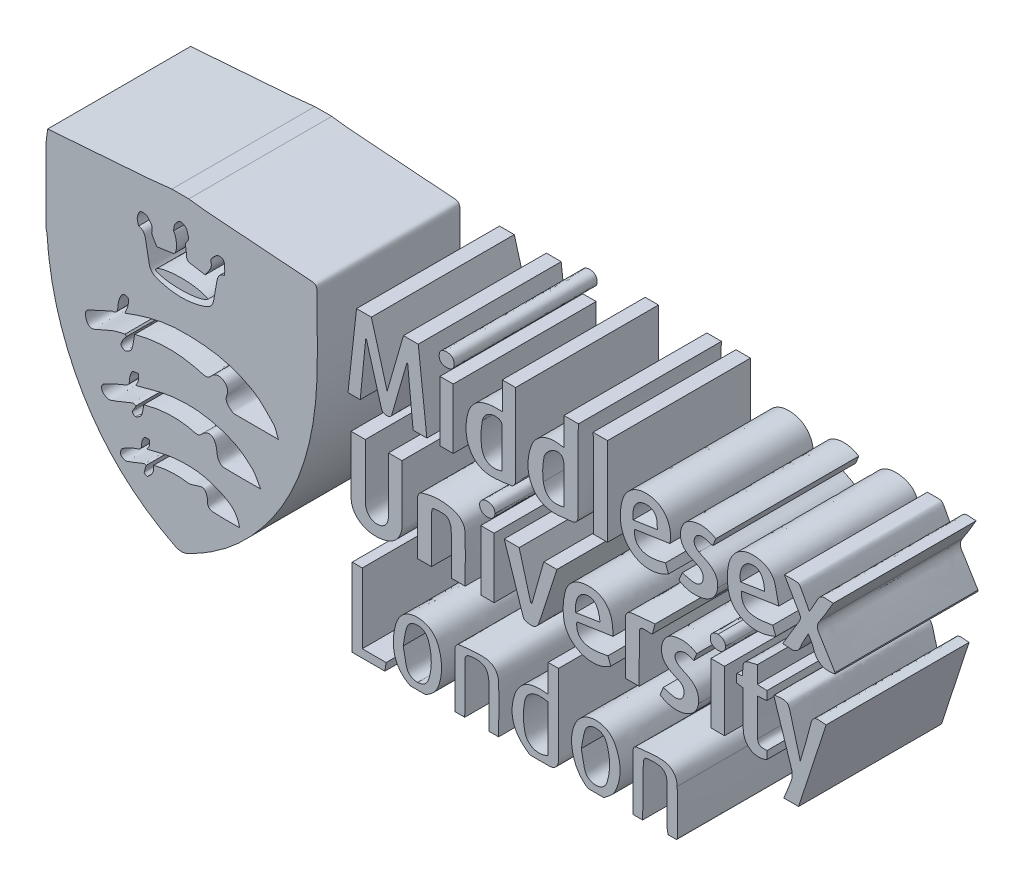
SolidWorks part; units mm, degrees
ref_plane "Front Plane" through (0, 0, 0) normal (0, 0, 1) x (1, 0, 0)
ref_plane "Top Plane" through (0, 0, 0) normal (0, 1, 0) x (1, 0, 0)
ref_plane "Right Plane" through (0, 0, 0) normal (1, 0, 0) x (0, 0, -1)
sketch "Model" plane through (0, 0, 0) normal (0, 0, 1) x (1, 0, 0)
  spline S0 degree 3 poles (174.4228, 110.9476) (174.5606, 110.6872) (174.6985, 110.5042) (174.7591, 110.2984) (174.9938, 109.5024) (175.5287, 109.2789) (176.2901, 109.4458) knots 92 92 92 92 93 93 93 94 94 94 94
  spline S1 degree 3 poles (173.8893, 109.9229) (174.0165, 110.2569) (174.2185, 110.5625) (174.4228, 110.9476) knots 91 91 91 91 92 92 92 92
  spline S2 degree 3 poles (172.6251, 109.454) (172.8108, 109.4445) (172.9346, 109.4503) (173.0539, 109.43) (173.4751, 109.3581) (173.7331, 109.5127) (173.8893, 109.9229) knots 89 89 89 89 90 90 90 91 91 91 91
  spline S3 degree 3 poles (173.7729, 111.368) (173.3875, 110.7517) (173.0235, 110.1221) (172.6251, 109.454) knots 88 88 88 88 89 89 89 89
  spline S4 degree 3 poles (172.7457, 113.6889) (173.1195, 113.0375) (173.4368, 112.4592) (173.7814, 111.8977) (173.9035, 111.6988) (173.8929, 111.5598) (173.7729, 111.368) knots 86 86 86 86 87 87 87 88 88 88 88
  spline S5 degree 3 poles (174.4932, 112.3338) (174.2779, 112.7438) (174.1029, 113.093) (173.9111, 113.4326) (173.855, 113.5319) (173.7581, 113.6671) (173.6677, 113.6773) (173.3856, 113.7091) (173.0976, 113.6889) (172.7457, 113.6889) knots 83 83 83 83 84 84 84 85 85 85 86 86 86 86
  spline S6 degree 3 poles (176.1595, 113.6612) (175.2657, 113.7417) (175.2671, 113.7409) (174.9095, 113.0736) (174.7857, 112.8426) (174.6527, 112.6165) (174.4932, 112.3338) knots 81 81 81 81 82 82 82 83 83 83 83
  spline S7 degree 3 poles (175.2088, 112.1108) (175.5437, 112.6021) (175.8336, 113.1241) (176.1595, 113.6612) knots 80 80 80 80 81 81 81 81
  spline S8 degree 3 poles (176.2901, 109.5304) (175.9311, 110.1153) (175.588, 110.7108) (175.2064, 111.2805) (175.006, 111.5798) (175.0052, 111.8119) (175.2088, 112.1108) knots 78 78 78 78 79 79 79 80 80 80 80
  spline S11 degree 3 poles (160.3728, 109.4654) (160.3728, 111.5413) (160.3728, 113.5839) (160.3728, 115.6264) knots 75 75 75 75 76 76 76 76
  spline S12 degree 3 poles (159.3992, 109.4654) (159.7501, 109.4654) (160.0504, 109.4654) (160.3728, 109.4654) knots 74 74 74 74 75 75 75 75
  spline S13 degree 3 poles (159.3568, 115.6264) (159.3709, 115.4595) (159.3971, 115.2926) (159.3974, 115.1257) (159.4004, 113.4059) (159.3992, 111.686) (159.3992, 109.9662) (159.3992, 109.8003) (159.3992, 109.6344) (159.3992, 109.4654) knots 71 71 71 71 72 72 72 73 73 73 74 74 74 74
  spline S15 degree 3 poles (154.8135, 111.5818) (154.7295, 110.4142) (155.3759, 109.4945) (156.3943, 109.3858) (156.8744, 109.3346) (157.3728, 109.4233) (157.8597, 109.4773) (158.1797, 109.5128) (158.3137, 109.6905) (158.3084, 110.0511) (158.285, 111.6437) (158.2964, 113.2368) (158.3002, 114.8297) (158.3009, 115.0953) (158.3266, 115.3609) (158.3408, 115.6264) knots 65 65 65 65 66 66 66 67 67 67 68 68 68 69 69 69 70 70 70 70
  spline S16 degree 3 poles (157.3248, 113.6773) (157.1356, 113.7017) (156.9969, 113.7232) (156.8576, 113.7368) (156.0697, 113.8138) (155.3479, 113.4198) (155.0538, 112.6876) (154.9149, 112.3417) (154.8404, 111.9554) (154.8135, 111.5818) knots 62 62 62 62 63 63 63 64 64 64 65 65 65 65
  spline S17 degree 3 poles (157.3248, 115.6264) (157.3248, 114.9831) (157.3248, 114.3399) (157.3248, 113.6773) knots 61 61 61 61 62 62 62 62
  spline S19 degree 3 poles (150.4908, 111.8155) (150.3546, 110.575) (150.8981, 109.5849) (151.921, 109.4274) (152.4861, 109.3404) (153.0888, 109.4634) (153.6687, 109.5374) (153.7772, 109.5513) (153.9386, 109.7813) (153.9395, 109.9125) (153.9527, 111.817) (153.9426, 113.7218) (153.9381, 115.6264) knots 56 56 56 56 57 57 57 58 58 58 59 59 59 60 60 60 60
  spline S20 degree 3 poles (153.0068, 113.7012) (151.3689, 113.7884) (150.6459, 113.2282) (150.4908, 111.8155) knots 55 55 55 55 56 56 56 56
  spline S21 degree 3 poles (153.0068, 115.6264) (153.0068, 114.9855) (153.0068, 114.3446) (153.0068, 113.7012) knots 54 54 54 54 55 55 55 55
  spline S23 degree 3 poles (121.0874, 108.8531) (121.1149, 108.7329) (121.1594, 108.6138) (121.1673, 108.4923) (121.2824, 106.7106) (121.6082, 104.9688) (122.2053, 103.2862) (123.6475, 99.2218) (126.1934, 96.1002) (130.0768, 94.1277) (130.4064, 93.9603) (130.6811, 93.9473) (131.0261, 94.114) (132.7644, 94.9538) (134.2736, 96.0965) (135.5682, 97.5178) (138.5327, 100.7727) (139.8486, 104.6871) (140.0355, 109.0137) (140.114, 110.8297) (140.0377, 112.6522) (140.0449, 114.4716) (140.0462, 114.7877) (139.9531, 114.9147) (139.6186, 114.9377) (137.2282, 115.102) (134.839, 115.2828) (132.45, 115.4663) (131.9913, 115.5016) (131.5353, 115.5722) (131.0781, 115.6264) knots 43 43 43 43 44 44 44 45 45 45 46 46 46 47 47 47 48 48 48 49 49 49 50 50 50 51 51 51 52 52 52 53 53 53 53
  spline S26 degree 3 poles (142.5081, 99.3333) (142.5081, 97.4962) (142.5081, 95.6817) (142.5081, 93.8671) knots 40 40 40 40 41 41 41 41
  spline S27 degree 3 poles (143.2124, 99.3333) (142.9542, 99.3333) (142.7483, 99.3333) (142.5081, 99.3333) knots 39 39 39 39 40 40 40 40
  spline S28 degree 3 poles (143.2124, 94.4354) (143.2124, 96.1023) (143.2124, 97.7159) (143.2124, 99.3333) knots 38 38 38 38 39 39 39 39
  spline S29 degree 3 poles (144.8804, 94.4354) (144.2895, 94.4354) (143.7758, 94.4354) (143.2124, 94.4354) knots 37 37 37 37 38 38 38 38
  spline S30 degree 3 poles (144.7941, 93.8671) (144.8197, 94.0356) (144.8453, 94.204) (144.8804, 94.4354) knots 36 36 36 36 37 37 37 37
  spline S32 degree 3 poles (147.5881, 93.8671) (148.0629, 94.0735) (148.4105, 94.4076) (148.5707, 94.9045) (148.8199, 95.6774) (148.8263, 96.4571) (148.555, 97.2258) (148.322, 97.8858) (147.8041, 98.2488) (147.1153, 98.2676) (146.4326, 98.2863) (145.887, 97.9454) (145.6323, 97.2937) (145.5211, 97.0091) (145.4516, 96.6999) (145.4155, 96.3957) (145.2709, 95.1793) (145.6611, 94.3457) (146.5721, 93.8671) knots 29 29 29 29 30 30 30 31 31 31 32 32 32 33 33 33 34 34 34 35 35 35 35
  spline S34 degree 3 poles (152.7528, 93.8671) (152.7585, 94.9489) (152.7868, 96.0313) (152.7612, 97.1123) (152.7469, 97.7142) (152.4166, 98.1234) (151.8172, 98.1738) (151.2005, 98.2257) (150.5684, 98.1294) (149.9474, 98.0591) (149.8501, 98.0481) (149.7038, 97.8319) (149.7025, 97.7092) (149.6889, 96.4287) (149.7003, 95.1478) (149.7048, 93.8671) knots 23 23 23 23 24 24 24 25 25 25 26 26 26 27 27 27 28 28 28 28
  spline S36 degree 3 poles (156.2142, 98.1705) (156.0514, 98.1828) (155.9393, 98.1894) (155.8277, 98.2001) (154.8095, 98.2973) (154.1122, 97.8257) (153.8313, 96.849) (153.4593, 95.5554) (153.8291, 94.5733) (154.9541, 93.8671) knots 19 19 19 19 20 20 20 21 21 21 22 22 22 22
  spline S37 degree 3 poles (156.2142, 100.1122) (156.2142, 99.4567) (156.2142, 98.8195) (156.2142, 98.1705) knots 18 18 18 18 19 19 19 19
  spline S38 degree 3 poles (156.9436, 100.1122) (156.6759, 100.1122) (156.47, 100.1122) (156.2142, 100.1122) knots 17 17 17 17 18 18 18 18
  spline S39 degree 3 poles (156.3934, 93.8671) (156.8995, 93.9891) (156.9648, 94.3302) (156.9557, 94.8027) (156.9244, 96.4217) (156.9436, 98.0417) (156.9436, 99.6613) (156.9436, 99.8102) (156.9436, 99.959) (156.9436, 100.1122) knots 14 14 14 14 15 15 15 16 16 16 17 17 17 17
  spline S41 degree 3 poles (160.1188, 93.8671) (160.3727, 94.0981) (160.7149, 94.2828) (160.8645, 94.5684) (161.3785, 95.5498) (161.3889, 96.5839) (160.8559, 97.5573) (160.3605, 98.4617) (158.9813, 98.5175) (158.3339, 97.7082) (157.4649, 96.6221) (157.8315, 94.5638) (159.0181, 93.8671) knots 9 9 9 9 10 10 10 11 11 11 12 12 12 13 13 13 13
  spline S43 degree 3 poles (165.2474, 97.1096) (165.2234, 97.7242) (164.8663, 98.13) (164.25, 98.1851) (163.6729, 98.2366) (163.0811, 98.1437) (162.4975, 98.0935) (162.2379, 98.0711) (162.1401, 97.9128) (162.1438, 97.6314) (162.1605, 96.3768) (162.1509, 95.1219) (162.1508, 93.8671) knots 4 4 4 4 5 5 5 6 6 6 7 7 7 8 8 8 8
  spline S44 degree 3 poles (165.1988, 93.8671) (165.2202, 93.9188) (165.2603, 93.9704) (165.2604, 94.0221) (165.2623, 95.0514) (165.2874, 96.0818) (165.2474, 97.1096) knots 2 2 2 2 3 3 3 4 4 4 4
  spline S47 degree 3 poles (143.0697, 109.457) (143.1991, 110.7616) (143.3262, 112.0442) (143.4533, 113.3268) knots 15 15 15 15 16 16 16 16
  spline S48 degree 3 poles (142.2133, 109.457) (142.5245, 109.457) (142.7844, 109.457) (143.0697, 109.457) knots 14 14 14 14 15 15 15 15
  spline S49 degree 3 poles (142.814, 114.8472) (142.6136, 113.049) (142.4146, 111.2634) (142.2133, 109.457) knots 13 13 13 13 14 14 14 14
  spline S50 degree 3 poles (143.8503, 114.8472) (143.4936, 114.8472) (143.1727, 114.8472) (142.814, 114.8472) knots 12 12 12 12 13 13 13 13
  spline S51 degree 3 poles (144.9531, 110.9127) (144.5616, 112.3095) (144.2055, 113.5799) (143.8503, 114.8472) knots 11 11 11 11 12 12 12 12
  spline S52 degree 3 poles (146.0946, 114.849) (145.7232, 113.5681) (145.3541, 112.2955) (144.9531, 110.9127) knots 10 10 10 10 11 11 11 11
  spline S53 degree 3 poles (147.1297, 114.849) (146.7576, 114.849) (146.4359, 114.849) (146.0946, 114.849) knots 9 9 9 9 10 10 10 10
  spline S54 degree 3 poles (147.7331, 109.4589) (147.5299, 111.274) (147.33, 113.0596) (147.1297, 114.849) knots 8 8 8 8 9 9 9 9
  spline S55 degree 3 poles (146.7711, 109.4589) (147.1034, 109.4589) (147.4055, 109.4589) (147.7331, 109.4589) knots 7 7 7 7 8 8 8 8
  spline S56 degree 3 poles (146.389, 113.3208) (146.5158, 112.0387) (146.6427, 110.7567) (146.7711, 109.4589) knots 6 6 6 6 7 7 7 7
  spline S57 degree 3 poles (146.3401, 113.3276) (146.3564, 113.3253) (146.3727, 113.323) (146.389, 113.3208) knots 5 5 5 5 6 6 6 6
  spline S58 degree 3 poles (143.5043, 113.3343) (143.8397, 112.1613) (144.1798, 110.9895) (144.5066, 109.8141) (144.5722, 109.5781) (144.6255, 109.4148) (144.9376, 109.4198) (145.2408, 109.4246) (145.2669, 109.6034) (145.3261, 109.8108) (145.6608, 110.984) (146.0015, 112.1555) (146.3401, 113.3276) knots 1 1 1 1 2 2 2 3 3 3 4 4 4 5 5 5 5
  spline S59 degree 3 poles (143.4533, 113.3268) (143.4703, 113.3293) (143.4873, 113.3318) (143.5043, 113.3343) knots 0 0 0 0 1 1 1 1
  spline S60 degree 3 poles (142.4263, 107.2195) (142.4263, 105.8316) (142.3913, 104.467) (142.4398, 103.1053) (142.4675, 102.3291) (143.1801, 101.7637) (144.0054, 101.7284) (145.0567, 101.6834) (145.78, 102.1367) (145.9626, 102.9567) (145.9778, 103.0251) (145.9877, 103.0963) (145.9878, 103.1662) (145.9893, 104.504) (145.9889, 105.8417) (145.9889, 107.2192) knots 9 9 9 9 10 10 10 11 11 11 12 12 12 13 13 13 14 14 14 14
  spline S61 degree 3 poles (143.4251, 107.2195) (143.0541, 107.2195) (142.7495, 107.2195) (142.4263, 107.2195) knots 8 8 8 8 9 9 9 9
  spline S62 degree 3 poles (145.0484, 107.2192) (145.0484, 107.0424) (145.0484, 106.8903) (145.0484, 106.7381) (145.0484, 105.611) (145.0544, 104.4838) (145.0455, 103.3567) (145.0415, 102.8558) (144.7347, 102.5276) (144.2885, 102.5056) (143.8277, 102.4829) (143.4842, 102.8064) (143.4391, 103.3131) (143.4255, 103.4671) (143.4259, 103.6226) (143.4257, 103.7775) (143.4246, 104.7778) (143.4251, 105.7782) (143.4251, 106.7785) (143.4251, 106.9268) (143.4251, 107.0752) (143.4251, 107.2195) knots 1 1 1 1 2 2 2 3 3 3 4 4 4 5 5 5 6 6 6 7 7 7 8 8 8 8
  spline S63 degree 3 poles (145.9889, 107.2192) (145.6549, 107.2192) (145.3677, 107.2192) (145.0484, 107.2192) knots 0 0 0 0 1 1 1 1
  spline S64 degree 3 poles (149.4511, 101.8273) (149.7999, 101.8273) (150.0796, 101.8273) (150.4118, 101.8273) knots 14 14 14 14 15 15 15 15
  spline S65 degree 3 poles (148.0536, 101.8302) (148.0536, 101.9991) (148.0536, 102.1508) (148.0536, 102.3025) (148.0537, 103.2181) (148.0497, 104.1337) (148.0585, 105.0492) (148.0598, 105.1786) (148.1119, 105.4139) (148.1602, 105.4192) (148.4731, 105.4535) (148.8179, 105.5113) (149.0979, 105.4105) (149.2663, 105.3499) (149.4256, 105.0205) (149.4352, 104.805) (149.4733, 103.9474) (149.451, 103.0872) (149.4511, 102.2279) (149.4511, 102.095) (149.4511, 101.9621) (149.4511, 101.8273) knots 7 7 7 7 8 8 8 9 9 9 10 10 10 11 11 11 12 12 12 13 13 13 14 14 14 14
  spline S66 degree 3 poles (147.0664, 101.8302) (147.419, 101.8302) (147.7107, 101.8302) (148.0536, 101.8302) knots 6 6 6 6 7 7 7 7
  spline S67 degree 3 poles (150.4118, 101.8273) (150.4118, 102.9392) (150.4381, 104.0084) (150.4009, 105.0753) (150.3819, 105.6177) (149.9908, 105.9274) (149.4873, 106.0538) (148.7588, 106.2368) (148.03, 106.173) (147.3255, 105.9353) (147.2082, 105.8957) (147.0813, 105.6789) (147.0779, 105.541) (147.0556, 104.6541) (147.0664, 103.7664) (147.0664, 102.879) (147.0664, 102.5326) (147.0664, 102.1863) (147.0664, 101.8302) knots 0 0 0 0 1 1 1 2 2 2 3 3 3 4 4 4 5 5 5 6 6 6 6
  spline S68 degree 3 poles (173.2553, 102.1372) (173.3156, 101.9425) (173.3027, 101.6941) (173.239, 101.4981) (173.0928, 101.0483) (172.8943, 100.6154) (172.7025, 100.1396) knots 10 10 10 10 11 11 11 12 12 12 12
  spline S69 degree 3 poles (172.1238, 105.6279) (172.5037, 104.4652) (172.8936, 103.3056) (173.2553, 102.1372) knots 9 9 9 9 10 10 10 10
  spline S70 degree 3 poles (172.0028, 106.0188) (172.0417, 105.8929) (172.0808, 105.7598) (172.1238, 105.6279) knots 8 8 8 8 9 9 9 9
  spline S71 degree 3 poles (173.8558, 102.9646) (173.6319, 103.8001) (173.4359, 104.529) (173.2413, 105.2583) (173.0009, 106.1593) (173.0015, 106.1595) (172.057, 106.0513) (172.0452, 106.05) (172.0346, 106.0383) (172.0028, 106.0188) knots 5 5 5 5 6 6 6 7 7 7 8 8 8 8
  spline S72 degree 3 poles (174.5794, 105.5349) (174.3932, 104.7054) (174.123, 103.8947) (173.8558, 102.9646) knots 4 4 4 4 5 5 5 5
  spline S73 degree 3 poles (175.6664, 106.0521) (175.5161, 106.0611) (175.4184, 106.0581) (175.3239, 106.0743) (174.8884, 106.1489) (174.6821, 105.9924) (174.5794, 105.5349) knots 2 2 2 2 3 3 3 4 4 4 4
  spline S74 degree 3 poles (173.7383, 100.1396) (174.3781, 102.1016) (175.0171, 104.0609) (175.6664, 106.0521) knots 1 1 1 1 2 2 2 2
  spline S75 degree 3 poles (172.7025, 100.1396) (173.0756, 100.1396) (173.3945, 100.1396) (173.7383, 100.1396) knots 0 0 0 0 1 1 1 1
  spline S76 degree 3 poles (162.2778, 111.206) (163.0927, 111.3276) (163.9122, 111.4499) (164.7298, 111.5719) knots 6 6 6 6 7 7 7 7
  spline S77 degree 3 poles (164.425, 110.2473) (162.9839, 109.8092) (162.142, 110.1883) (162.2778, 111.206) knots 5 5 5 5 6 6 6 6
  spline S78 degree 3 poles (164.6399, 109.6805) (164.5693, 109.8665) (164.4967, 110.058) (164.425, 110.2473) knots 4 4 4 4 5 5 5 5
  spline S79 degree 3 poles (164.7298, 111.5719) (164.9553, 112.5531) (164.4514, 113.4964) (163.5874, 113.7173) (162.5646, 113.9789) (161.6632, 113.4866) (161.3887, 112.4766) (161.2944, 112.1297) (161.2574, 111.7535) (161.2703, 111.3934) (161.3345, 109.6077) (163.0603, 108.7212) (164.6399, 109.6805) knots 0 0 0 0 1 1 1 2 2 2 3 3 3 4 4 4 4
  spline S80 degree 3 poles (169.7327, 111.2022) (170.5641, 111.3258) (171.399, 111.4499) (172.3562, 111.5922) knots 8 8 8 8 9 9 9 9
  spline S81 degree 3 poles (171.9257, 110.2205) (170.2967, 109.9082) (169.716, 110.1672) (169.7327, 111.2022) knots 7 7 7 7 8 8 8 8
  spline S82 degree 3 poles (172.1459, 109.6451) (172.0623, 109.8636) (171.9931, 110.0444) (171.9257, 110.2205) knots 6 6 6 6 7 7 7 7
  spline S83 degree 3 poles (169.7348, 109.5758) (170.5307, 109.1814) (171.3373, 109.2981) (172.1459, 109.6451) knots 5 5 5 5 6 6 6 6
  spline S84 degree 3 poles (168.8439, 112.3798) (168.7731, 112.068) (168.754, 111.7377) (168.7592, 111.4167) (168.7717, 110.6436) (168.9919, 109.944) (169.7348, 109.5758) knots 3 3 3 3 4 4 4 5 5 5 5
  spline S85 degree 3 poles (172.3562, 111.5922) (172.2528, 112.0546) (172.1953, 112.4854) (172.0561, 112.888) (171.8987, 113.3432) (171.5315, 113.605) (171.0617, 113.721) (170.0011, 113.983) (169.0851, 113.4419) (168.8439, 112.3798) knots 0 0 0 0 1 1 1 2 2 2 3 3 3 3
  spline S86 degree 3 poles (158.2238, 103.5789) (159.0527, 103.7026) (159.8851, 103.8269) (160.7585, 103.9573) knots 7 7 7 7 8 8 8 8
  spline S87 degree 3 poles (160.4004, 102.6055) (158.8527, 102.239) (158.1293, 102.5675) (158.2238, 103.5789) knots 6 6 6 6 7 7 7 7
  spline S88 degree 3 poles (160.5977, 102.0737) (160.5318, 102.2512) (160.4651, 102.4311) (160.4004, 102.6055) knots 5 5 5 5 6 6 6 6
  spline S89 degree 3 poles (157.4007, 104.973) (157.2609, 104.4179) (157.2153, 103.7912) (157.319, 103.2321) (157.5828, 101.8093) (159.4073, 101.1891) (160.5977, 102.0737) knots 3 3 3 3 4 4 4 5 5 5 5
  spline S90 degree 3 poles (160.7585, 103.9573) (160.7436, 104.2014) (160.7419, 104.4243) (160.7144, 104.644) (160.6053, 105.5151) (160.0872, 106.0604) (159.3059, 106.1385) (158.3658, 106.2325) (157.6173, 105.8321) (157.4007, 104.973) knots 0 0 0 0 1 1 1 2 2 2 3 3 3 3
  spline S91 degree 3 poles (154.1902, 106.0545) (153.8491, 106.0545) (153.5289, 106.0545) (153.1442, 106.0545) knots 9 9 9 9 10 10 10 10
  spline S92 degree 3 poles (154.9966, 103.1258) (154.7288, 104.0982) (154.4611, 105.0706) (154.1902, 106.0545) knots 8 8 8 8 9 9 9 9
  spline S93 degree 3 poles (155.0817, 103.1146) (155.0533, 103.1184) (155.0249, 103.1221) (154.9966, 103.1258) knots 7 7 7 7 8 8 8 8
  spline S94 degree 3 poles (155.9096, 106.0499) (155.6301, 105.0587) (155.3559, 104.0867) (155.0817, 103.1146) knots 6 6 6 6 7 7 7 7
  spline S95 degree 3 poles (156.8286, 106.0499) (156.4967, 106.0499) (156.2066, 106.0499) (155.9096, 106.0499) knots 5 5 5 5 6 6 6 6
  spline S96 degree 3 poles (153.1442, 106.0545) (153.5967, 104.6615) (154.0285, 103.3249) (154.4702, 101.9916) (154.4944, 101.9186) (154.5937, 101.8386) (154.6716, 101.8205) (155.2588, 101.6842) (155.4678, 101.8086) (155.6465, 102.3757) (155.6803, 102.483) (155.7199, 102.5885) (155.7542, 102.6956) (156.1099, 103.8049) (156.465, 104.9144) (156.8286, 106.0499) knots 0 0 0 0 1 1 1 2 2 2 3 3 3 4 4 4 5 5 5 5
  spline S97 degree 3 poles (169.4122, 105.4641) (169.5644, 105.4359) (169.6979, 105.4112) (169.8588, 105.3814) knots 13 13 13 13 14 14 14 14
  spline S98 degree 3 poles (169.4122, 106.0377) (169.4122, 105.8338) (169.4122, 105.6559) (169.4122, 105.4641) knots 12 12 12 12 13 13 13 13
  spline S99 degree 3 poles (169.8136, 106.0988) (169.6833, 106.079) (169.5507, 106.0588) (169.4122, 106.0377) knots 11 11 11 11 12 12 12 12
  spline S100 degree 3 poles (170.8518, 107.2904) (170.5087, 107.1863) (170.1208, 107.1806) (169.953, 106.9856) (169.7898, 106.7958) (169.8521, 106.4121) (169.8136, 106.0988) knots 9 9 9 9 10 10 10 11 11 11 11
  spline S101 degree 3 poles (170.8518, 106.0966) (170.8518, 106.4956) (170.8518, 106.8574) (170.8518, 107.2904) knots 8 8 8 8 9 9 9 9
  spline S102 degree 3 poles (171.523, 106.0561) (171.2944, 106.0699) (171.09, 106.0822) (170.8518, 106.0966) knots 7 7 7 7 8 8 8 8
  spline S103 degree 3 poles (171.523, 105.4526) (171.523, 105.6622) (171.523, 105.8524) (171.523, 106.0561) knots 6 6 6 6 7 7 7 7
  spline S104 degree 3 poles (170.8669, 105.3939) (171.1062, 105.4153) (171.3122, 105.4338) (171.523, 105.4526) knots 5 5 5 5 6 6 6 6
  spline S105 degree 3 poles (170.8753, 102.8085) (170.8487, 103.6647) (170.8669, 104.5222) (170.8669, 105.3939) knots 4 4 4 4 5 5 5 5
  spline S106 degree 3 poles (171.5262, 102.4241) (171.2039, 102.4049) (170.887, 102.4302) (170.8753, 102.8085) knots 3 3 3 3 4 4 4 4
  spline S107 degree 3 poles (171.5262, 101.88) (171.5262, 102.0608) (171.5262, 102.2397) (171.5262, 102.4241) knots 2 2 2 2 3 3 3 3
  spline S108 degree 3 poles (169.8588, 105.3814) (169.8588, 104.5392) (169.8373, 103.7078) (169.8646, 102.8779) (169.895, 101.9531) (170.6885, 101.4922) (171.5262, 101.88) knots 0 0 0 0 1 1 1 2 2 2 2
  spline S109 degree 3 poles (165.6032, 110.2396) (165.5276, 110.06) (165.4521, 109.8803) (165.3626, 109.6675) knots 15 15 15 15 16 16 16 16
  spline S110 degree 3 poles (167.038, 110.4709) (166.9416, 110.1377) (166.6583, 110.0221) (166.3373, 110.0594) (166.0948, 110.0876) (165.8591, 110.1745) (165.6032, 110.2396) knots 13 13 13 13 14 14 14 15 15 15 15
  spline S111 degree 3 poles (167.9458, 113.4697) (167.4333, 113.7859) (166.9148, 113.8507) (166.3787, 113.706) (165.8498, 113.5634) (165.5522, 113.192) (165.4775, 112.6509) (165.4108, 112.1677) (165.6524, 111.7384) (166.1352, 111.479) (166.3082, 111.3861) (166.4927, 111.3146) (166.6711, 111.2314) (167, 111.0779) (167.1364, 110.8108) (167.038, 110.4709) knots 8 8 8 8 9 9 9 10 10 10 11 11 11 12 12 12 13 13 13 13
  spline S112 degree 3 poles (167.7359, 112.9407) (167.8082, 113.1231) (167.8739, 113.2886) (167.9458, 113.4697) knots 7 7 7 7 8 8 8 8
  spline S113 degree 3 poles (166.7625, 112.0718) (166.4847, 112.2308) (166.3593, 112.4702) (166.4785, 112.7822) (166.5921, 113.0795) (166.8482, 113.158) (167.1352, 113.1116) (167.3347, 113.0793) (167.5269, 113.0019) (167.7359, 112.9407) knots 4 4 4 4 5 5 5 6 6 6 7 7 7 7
  spline S114 degree 3 poles (168.0745, 110.5419) (168.129, 111.126) (167.8713, 111.5327) (167.2554, 111.8326) (167.0912, 111.9126) (166.9206, 111.9813) (166.7625, 112.0718) knots 2 2 2 2 3 3 3 4 4 4 4
  spline S115 degree 3 poles (165.3626, 109.6675) (165.8952, 109.3428) (166.4362, 109.293) (166.9865, 109.4028) (167.6068, 109.5266) (168.0226, 109.9862) (168.0745, 110.5419) knots 0 0 0 0 1 1 1 2 2 2 2
  spline S116 degree 3 poles (164.1649, 105.0812) (164.0841, 104.5257) (164.2959, 104.121) (164.8269, 103.8385) (165, 103.7464) (165.185, 103.6769) (165.3626, 103.5931) (165.6792, 103.4438) (165.7844, 103.1795) (165.7031, 102.8592) (165.6163, 102.5168) (165.3379, 102.399) (165.0189, 102.4323) (164.7751, 102.4577) (164.5384, 102.5516) (164.2712, 102.6223) knots 11 11 11 11 12 12 12 13 13 13 14 14 14 15 15 15 16 16 16 16
  spline S117 degree 3 poles (166.6082, 105.835) (166.1466, 106.1573) (165.6485, 106.2036) (165.1412, 106.1101) (164.5984, 106.01) (164.2415, 105.6078) (164.1649, 105.0812) knots 9 9 9 9 10 10 10 11 11 11 11
  spline S118 degree 3 poles (166.4054, 105.3173) (166.4725, 105.4885) (166.5381, 105.6562) (166.6082, 105.835) knots 8 8 8 8 9 9 9 9
  spline S119 degree 3 poles (165.1512, 105.1356) (165.2623, 105.3127) (165.5326, 105.4483) (165.7507, 105.4828) (165.9481, 105.514) (166.1711, 105.383) (166.4054, 105.3173) knots 6 6 6 6 7 7 7 8 8 8 8
  spline S120 degree 3 poles (166.7298, 102.8627) (166.7985, 103.4768) (166.5676, 103.884) (165.9734, 104.187) (165.7858, 104.2826) (165.5851, 104.3549) (165.4051, 104.4626) (165.1482, 104.6163) (164.9909, 104.88) (165.1512, 105.1356) knots 3 3 3 3 4 4 4 5 5 5 6 6 6 6
  spline S121 degree 3 poles (164.0491, 102.0627) (164.5345, 101.738) (165.1883, 101.6376) (165.7271, 101.7918) (166.2998, 101.9558) (166.673, 102.3543) (166.7298, 102.8627) knots 1 1 1 1 2 2 2 3 3 3 3
  spline S122 degree 3 poles (164.2712, 102.6223) (164.1987, 102.4397) (164.1227, 102.2482) (164.0491, 102.0627) knots 0 0 0 0 1 1 1 1
  spline S123 degree 3 poles (163.5049, 105.4831) (163.5584, 105.6747) (163.6145, 105.8756) (163.7008, 106.1847) knots 8 8 8 8 9 9 9 9
  spline S124 degree 3 poles (162.5878, 101.8487) (162.5878, 102.8275) (162.5879, 103.7697) (162.5878, 104.712) (162.5877, 105.5188) (162.5877, 105.5185) (163.4082, 105.4546) (163.4336, 105.4526) (163.4605, 105.4695) (163.5049, 105.4831) knots 5 5 5 5 6 6 6 7 7 7 8 8 8 8
  spline S125 degree 3 poles (161.629, 101.8487) (161.9756, 101.8487) (162.2728, 101.8487) (162.5878, 101.8487) knots 4 4 4 4 5 5 5 5
  spline S126 degree 3 poles (163.7008, 106.1847) (163.1455, 106.1325) (162.6577, 106.0938) (162.1717, 106.0388) (161.7643, 105.9928) (161.568, 105.794) (161.6194, 105.3434) (161.6653, 104.9406) (161.629, 104.5284) (161.629, 104.1203) (161.629, 103.3647) (161.629, 102.6092) (161.629, 101.8487) knots 0 0 0 0 1 1 1 2 2 2 3 3 3 4 4 4 4
  spline S127 degree 3 poles (148.6468, 109.4497) (148.9663, 109.4497) (149.2575, 109.4497) (149.5774, 109.4497) knots 3 3 3 3 4 4 4 4
  spline S128 degree 3 poles (148.6468, 113.6587) (148.6468, 112.2386) (148.6468, 110.8528) (148.6468, 109.4497) knots 2 2 2 2 3 3 3 3
  spline S129 degree 3 poles (149.5774, 113.6587) (149.2485, 113.6587) (148.9484, 113.6587) (148.6468, 113.6587) knots 1 1 1 1 2 2 2 2
  spline S130 degree 3 poles (149.5774, 109.4497) (149.5774, 110.8863) (149.5774, 112.2721) (149.5774, 113.6587) knots 0 0 0 0 1 1 1 1
  spline S131 degree 3 poles (152.434, 101.8356) (152.434, 103.2477) (152.434, 104.6363) (152.434, 106.048) knots 3 3 3 3 4 4 4 4
  spline S132 degree 3 poles (151.504, 101.8356) (151.8306, 101.8356) (152.1216, 101.8356) (152.434, 101.8356) knots 2 2 2 2 3 3 3 3
  spline S133 degree 3 poles (151.504, 106.048) (151.504, 104.6256) (151.504, 103.2283) (151.504, 101.8356) knots 1 1 1 1 2 2 2 2
  spline S134 degree 3 poles (152.434, 106.048) (152.1112, 106.048) (151.8106, 106.048) (151.504, 106.048) knots 0 0 0 0 1 1 1 1
  spline S135 degree 3 poles (167.6062, 101.8374) (167.9305, 101.8374) (168.2327, 101.8374) (168.5596, 101.8374) knots 3 3 3 3 4 4 4 4
  spline S136 degree 3 poles (167.6062, 106.0469) (167.6062, 104.6348) (167.6062, 103.2488) (167.6062, 101.8374) knots 2 2 2 2 3 3 3 3
  spline S137 degree 3 poles (168.5596, 106.0469) (168.2314, 106.0469) (167.9293, 106.0469) (167.6062, 106.0469) knots 1 1 1 1 2 2 2 2
  spline S138 degree 3 poles (168.5596, 101.8374) (168.5596, 103.2659) (168.5596, 104.6531) (168.5596, 106.0469) knots 0 0 0 0 1 1 1 1
  spline S139 degree 3 poles (168.622, 107.2818) (168.6011, 107.6075) (168.3907, 107.7343) (168.0953, 107.756) knots 3 3 3 3 4 4 4 4
  spline S140 degree 3 poles (168.0953, 107.756) (167.7865, 107.7364) (167.5737, 107.6018) (167.5638, 107.2788) (167.5536, 106.9473) (167.7769, 106.8098) (168.0725, 106.7884) (168.3901, 106.7653) (168.6403, 106.9944) (168.622, 107.2818) knots 0 0 0 0 1 1 1 2 2 2 3 3 3 3
  spline S141 degree 3 poles (151.4225, 107.2675) (151.4435, 106.95) (151.6536, 106.8098) (151.9548, 106.7858) knots 3 3 3 3 4 4 4 4
  spline S142 degree 3 poles (152.4938, 107.2553) (152.4907, 107.579) (152.2943, 107.7307) (151.9881, 107.7499) (151.6723, 107.7698) (151.4038, 107.5494) (151.4225, 107.2675) knots 1 1 1 1 2 2 2 3 3 3 3
  spline S143 degree 3 poles (151.9548, 106.7858) (152.2495, 106.782) (152.4963, 106.9864) (152.4938, 107.2553) knots 0 0 0 0 1 1 1 1
  spline S144 degree 3 poles (148.5943, 114.8873) (148.5961, 114.5435) (148.8248, 114.4354) (149.0984, 114.4173) knots 3 3 3 3 4 4 4 4
  spline S145 degree 3 poles (149.0984, 114.4173) (149.4384, 114.4325) (149.6504, 114.5822) (149.6439, 114.9061) (149.6374, 115.229) (149.4156, 115.3817) (149.1072, 115.376) (148.8001, 115.3703) (148.5926, 115.2208) (148.5943, 114.8873) knots 0 0 0 0 1 1 1 2 2 2 3 3 3 3
  spline S146 degree 3 poles (129.8928, 115.6264) (130.2879, 115.6264) (130.683, 115.6264) (131.0781, 115.6264) knots 14 14 14 14 15 15 15 15
  spline S147 degree 3 poles (121.2054, 114.9269) (123.5616, 115.1023) (125.8936, 115.2726) (128.225, 115.4519) (128.7821, 115.4948) (129.3369, 115.5675) (129.8928, 115.6264) knots 12 12 12 12 13 13 13 14 14 14 14
  spline S148 degree 3 poles (121.0874, 114.0178) (121.1262, 114.3162) (121.1649, 114.6147) (121.2054, 114.9269) knots 11 11 11 11 12 12 12 12
  spline S149 degree 3 poles (121.0874, 108.8531) (121.0874, 110.5747) (121.0874, 112.2962) (121.0874, 114.0178) knots 10 10 10 10 11 11 11 11
  spline S150 degree 3 poles (131.0781, 115.6264) (131.5353, 115.5722) (131.9913, 115.5016) (132.45, 115.4663) (134.839, 115.2828) (137.2282, 115.102) (139.6186, 114.9377) (139.9531, 114.9147) (140.0462, 114.7877) (140.0449, 114.4716) (140.0377, 112.6522) (140.114, 110.8297) (140.0355, 109.0137) (139.8486, 104.6871) (138.5327, 100.7727) (135.5682, 97.5178) (134.2736, 96.0965) (132.7644, 94.9538) (131.0261, 94.114) (130.6811, 93.9473) (130.4064, 93.9603) (130.0768, 94.1277) (126.1934, 96.1002) (123.6475, 99.2218) (122.2053, 103.2862) (121.6082, 104.9688) (121.2824, 106.7106) (121.1673, 108.4923) (121.1594, 108.6138) (121.1149, 108.7329) (121.0874, 108.8531) knots 0 0 0 0 1 1 1 2 2 2 3 3 3 4 4 4 5 5 5 6 6 6 7 7 7 8 8 8 9 9 9 10 10 10 10
  spline S151 degree 3 poles (137.3453, 104.1863) (137.2131, 104.493) (137.1687, 104.77) (137.0087, 104.9347) (136.5526, 105.4043) (136.1058, 105.9224) (135.5541, 106.252) (134.0194, 107.1689) (132.2958, 107.3764) (130.5418, 107.3499) (129.2168, 107.3299) (127.9554, 106.9787) (126.6028, 106.4676) knots 24 24 24 24 25 25 25 26 26 26 27 27 27 28 28 28 28
  spline S152 degree 3 poles (127.2904, 105.5254) (128.7915, 105.9259) (130.3735, 105.9899) (131.9546, 105.5246) (132.2362, 105.4418) (132.4318, 105.4148) (132.6451, 105.6712) (132.8406, 105.9062) (133.1338, 106.0335) (133.4426, 105.871) (133.765, 105.7013) (133.8595, 105.3671) (133.7444, 105.0698) (133.5832, 104.6536) (133.8242, 104.4728) (134.0751, 104.2671) (134.1256, 104.2257) (134.1992, 104.19) (134.2623, 104.1897) (135.2577, 104.1849) (136.2531, 104.1863) (137.3453, 104.1863) knots 17 17 17 17 18 18 18 19 19 19 20 20 20 21 21 21 22 22 22 23 23 23 24 24 24 24
  spline S153 degree 3 poles (126.716, 105.0975) (126.6294, 104.9873) (126.5278, 104.8853) (126.4605, 104.7643) (126.3981, 104.6521) (126.3136, 104.4992) (126.3472, 104.4015) (126.3802, 104.3056) (126.5719, 104.1798) (126.6545, 104.2036) (126.8144, 104.2497) (127.0236, 104.3632) (127.0745, 104.5) (127.1876, 104.8039) (127.2155, 105.1394) (127.2904, 105.5254) knots 12 12 12 12 13 13 13 14 14 14 15 15 15 16 16 16 17 17 17 17
  spline S154 degree 3 poles (126.6265, 105.2109) (126.6564, 105.1731) (126.6862, 105.1353) (126.716, 105.0975) knots 11 11 11 11 12 12 12 12
  spline S155 degree 3 poles (126.6028, 106.4676) (126.6973, 106.6942) (126.773, 106.8253) (126.8053, 106.9663) (126.8432, 107.1319) (126.9213, 107.3718) (126.8442, 107.463) (126.6733, 107.6654) (126.4232, 107.5673) (126.3195, 107.3634) (126.2036, 107.1354) (126.131, 106.8663) (126.1169, 106.6108) (126.1025, 106.3494) (126.0583, 106.1793) (125.7668, 106.1523) (125.6879, 106.145) (125.6111, 106.1006) (125.5363, 106.0667) (125.0689, 105.8546) (124.6084, 105.6258) (124.1335, 105.4321) (123.7856, 105.2903) (123.8133, 105.0238) (123.891, 104.7664) (123.9701, 104.5043) (124.1681, 104.308) (124.4678, 104.4212) (124.9063, 104.5868) (125.3222, 104.8122) (125.7599, 104.9804) (126.0373, 105.087) (126.3369, 105.1361) (126.6265, 105.2109) knots 0 0 0 0 1 1 1 2 2 2 3 3 3 4 4 4 5 5 5 6 6 6 7 7 7 8 8 8 9 9 9 10 10 10 11 11 11 11
  spline S156 degree 3 poles (127.3962, 101.2522) (127.3673, 101.185) (127.3592, 101.1579) (127.3449, 101.1345) (127.2655, 101.0039) (127.1657, 100.8806) (127.1181, 100.7395) (127.1069, 100.7064) (127.3003, 100.5427) (127.3481, 100.5626) (127.5047, 100.6278) (127.6983, 100.7202) (127.7655, 100.8572) (127.8659, 101.0615) (127.8709, 101.3128) (127.9241, 101.5826) knots 20 20 20 20 21 21 21 22 22 22 23 23 23 24 24 24 25 25 25 25
  spline S157 degree 3 poles (127.5432, 103.2824) (127.396, 103.2492) (127.1821, 103.2639) (127.1164, 103.1722) (127.0026, 103.0135) (126.9396, 102.7908) (126.9307, 102.5916) (126.92, 102.352) (126.8751, 102.2209) (126.6214, 102.1257) (126.1304, 101.9412) (125.6552, 101.7095) (125.1877, 101.4697) (124.9392, 101.3423) (124.9171, 101.079) (125.0773, 100.8919) (125.1862, 100.7648) (125.4446, 100.642) (125.5828, 100.6858) (126.1126, 100.8534) (126.6191, 101.0938) (127.1394, 101.2939) (127.2067, 101.3198) (127.3035, 101.2692) (127.3962, 101.2522) knots 12 12 12 12 13 13 13 14 14 14 15 15 15 16 16 16 17 17 17 18 18 18 19 19 19 20 20 20 20
  spline S158 degree 3 poles (127.36, 102.4627) (127.4543, 102.648) (127.5324, 102.7438) (127.5496, 102.8494) (127.5723, 102.9897) (127.5476, 103.1377) (127.5432, 103.2824) knots 10 10 10 10 11 11 11 12 12 12 12
  spline S159 degree 3 poles (136.1044, 100.5602) (135.8679, 100.9509) (135.748, 101.2844) (135.5175, 101.4993) (135.1414, 101.8499) (134.7293, 102.2007) (134.2689, 102.4148) (132.7173, 103.1365) (131.0772, 103.3005) (129.3995, 102.9776) (128.7466, 102.8519) (128.1076, 102.6539) (127.36, 102.4627) knots 6 6 6 6 7 7 7 8 8 8 9 9 9 10 10 10 10
  spline S160 degree 3 poles (127.9241, 101.5826) (129.069, 101.8871) (130.2457, 102.0167) (131.4354, 101.6877) (131.6662, 101.6239) (131.8183, 101.6354) (131.9867, 101.8283) (132.1935, 102.0652) (132.5185, 102.2154) (132.7703, 101.9975) (132.9447, 101.8465) (133.026, 101.5231) (133.0416, 101.2701) (133.0607, 100.9595) (133.2258, 100.5822) (133.5342, 100.5705) (134.3424, 100.5399) (135.1525, 100.5602) (136.1044, 100.5602) knots 0 0 0 0 1 1 1 2 2 2 3 3 3 4 4 4 5 5 5 6 6 6 6
  spline S161 degree 3 poles (127.5652, 112.2242) (127.9289, 112.1774) (128.0194, 111.8876) (128.0756, 111.5682) (128.1416, 111.1938) (128.2278, 110.8223) (128.2767, 110.4458) (128.3254, 110.0697) (128.5101, 109.8154) (128.8625, 109.6916) (129.9927, 109.2947) (131.1269, 109.2958) (132.2568, 109.6892) (132.5873, 109.8043) (132.7822, 110.0366) (132.8276, 110.4038) (132.876, 110.7944) (132.967, 111.1796) (133.0333, 111.5681) (133.0883, 111.8905) (133.1852, 112.1748) (133.5654, 112.223) knots 20 20 20 20 21 21 21 22 22 22 23 23 23 24 24 24 25 25 25 26 26 26 27 27 27 27
  spline S162 degree 3 poles (128.8423, 111.6071) (128.7152, 111.8658) (128.4347, 112.1688) (128.493, 112.3771) (128.5969, 112.7486) (128.3534, 112.8976) (128.2038, 113.0812) (128.1179, 113.1865) (127.8218, 113.2301) (127.6955, 113.162) (127.569, 113.0939) (127.5013, 112.858) (127.4729, 112.6849) (127.4505, 112.5483) (127.527, 112.3955) (127.5652, 112.2242) knots 15 15 15 15 16 16 16 17 17 17 18 18 18 19 19 19 20 20 20 20
  spline S163 degree 3 poles (130.0066, 113.1504) (130.2363, 112.8776) (130.2976, 112.1016) (130.1, 111.8497) (130.0629, 111.8023) (129.984, 111.774) (129.92, 111.7638) (129.5768, 111.709) (129.2322, 111.6628) (128.8423, 111.6071) knots 12 12 12 12 13 13 13 14 14 14 15 15 15 15
  spline S164 degree 3 poles (132.2245, 111.5936) (131.9601, 111.6435) (131.7149, 111.703) (131.4661, 111.733) (131.2008, 111.7651) (130.9091, 111.7248) (130.9143, 112.1342) (130.9177, 112.3962) (130.7756, 112.7655) (130.9, 112.8988) (131.1646, 113.1822) (131.0169, 113.4318) (130.9474, 113.662) (130.906, 113.7995) (130.6612, 113.9653) (130.5172, 113.957) (130.374, 113.9488) (130.2108, 113.7588) (130.1155, 113.6105) (130.0352, 113.4854) (130.0396, 113.3058) (130.0066, 113.1504) knots 5 5 5 5 6 6 6 7 7 7 8 8 8 9 9 9 10 10 10 11 11 11 12 12 12 12
  spline S165 degree 3 poles (133.5654, 112.223) (133.5774, 112.3475) (133.6027, 112.4539) (133.5943, 112.5577) (133.5786, 112.7509) (133.5927, 112.9741) (133.4975, 113.1228) (133.4414, 113.2102) (133.1458, 113.2522) (133.0515, 113.1844) (132.8629, 113.049) (132.5762, 112.7724) (132.6166, 112.645) (132.7736, 112.1503) (132.3877, 111.9334) (132.2245, 111.5936) knots 0 0 0 0 1 1 1 2 2 2 3 3 3 4 4 4 5 5 5 5
  spline S166 degree 3 poles (128.6151, 98.2506) (129.403, 98.4603) (130.2043, 98.5239) (131.0251, 98.3853) (131.1767, 98.3597) (131.3478, 98.4488) (131.5097, 98.4859) (131.7157, 98.5331) (131.9848, 98.6825) (132.1112, 98.6033) (132.2686, 98.5048) (132.398, 98.2092) (132.379, 98.0144) (132.3444, 97.6599) (132.5497, 97.5132) (132.7885, 97.4965) (133.3883, 97.4547) (133.9929, 97.4827) (134.6262, 97.4827) knots 17 17 17 17 18 18 18 19 19 19 20 20 20 21 21 21 22 22 22 23 23 23 23
  spline S167 degree 3 poles (128.0969, 97.9939) (128.0393, 97.7986) (127.9779, 97.6409) (127.9574, 97.4781) (127.9535, 97.4464) (128.1553, 97.3389) (128.1825, 97.3616) (128.3246, 97.4804) (128.4722, 97.6135) (128.5562, 97.7739) (128.6217, 97.8989) (128.5969, 98.0712) (128.6151, 98.2506) knots 13 13 13 13 14 14 14 15 15 15 16 16 16 17 17 17 17
  spline S168 degree 3 poles (128.3062, 99.6781) (128.1807, 99.6534) (127.9973, 99.6707) (127.9423, 99.5949) (127.8427, 99.4576) (127.7793, 99.2658) (127.7747, 99.0948) (127.7685, 98.8679) (127.7308, 98.7584) (127.4791, 98.6821) (127.1167, 98.5721) (126.7677, 98.392) (126.4454, 98.1902) (126.3419, 98.1254) (126.2663, 97.8652) (126.3144, 97.7527) (126.3609, 97.6438) (126.6085, 97.524) (126.7232, 97.5583) (127.1406, 97.683) (127.5377, 97.8746) (127.9471, 98.0287) (128.001, 98.049) (128.0817, 97.9979) (128.0969, 97.9939) knots 5 5 5 5 6 6 6 7 7 7 8 8 8 9 9 9 10 10 10 11 11 11 12 12 12 13 13 13 13
  spline S169 degree 3 poles (128.1494, 99.003) (128.2297, 99.1378) (128.3082, 99.2176) (128.3235, 99.3082) (128.3438, 99.4271) (128.3143, 99.5544) (128.3062, 99.6781) knots 3 3 3 3 4 4 4 5 5 5 5
  spline S170 degree 3 poles (134.6262, 97.4827) (134.5029, 98.0939) (134.2271, 98.4626) (133.6197, 98.7938) (132.5057, 99.4012) (131.2962, 99.5479) (130.0583, 99.4102) (129.4421, 99.3417) (128.839, 99.1543) (128.1494, 99.003) knots 0 0 0 0 1 1 1 2 2 2 3 3 3 3
  spline S171 degree 3 poles (157.3248, 115.6264) (157.6634, 115.6264) (158.0021, 115.6264) (158.3408, 115.6264) knots 9 9 9 9 10 10 10 10
  spline S172 degree 3 poles (157.3248, 113.6773) (157.3248, 114.3399) (157.3248, 114.9831) (157.3248, 115.6264) knots 8 8 8 8 9 9 9 9
  spline S173 degree 3 poles (154.8135, 111.5818) (154.8404, 111.9554) (154.9149, 112.3417) (155.0538, 112.6876) (155.3479, 113.4198) (156.0697, 113.8138) (156.8576, 113.7368) (156.9969, 113.7232) (157.1356, 113.7017) (157.3248, 113.6773) knots 5 5 5 5 6 6 6 7 7 7 8 8 8 8
  spline S174 degree 3 poles (158.3408, 115.6264) (158.3266, 115.3609) (158.3009, 115.0953) (158.3002, 114.8297) (158.2964, 113.2368) (158.285, 111.6437) (158.3084, 110.0511) (158.3137, 109.6905) (158.1797, 109.5128) (157.8597, 109.4773) (157.3728, 109.4233) (156.8744, 109.3346) (156.3943, 109.3858) (155.3759, 109.4945) (154.7295, 110.4142) (154.8135, 111.5818) knots 0 0 0 0 1 1 1 2 2 2 3 3 3 4 4 4 5 5 5 5
  spline S175 degree 3 poles (155.8802, 110.8882) (156.0038, 110.1074) (156.5093, 109.8459) (157.3251, 110.0795) knots 4 4 4 4 5 5 5 5
  spline S176 degree 3 poles (157.3251, 110.0795) (157.3251, 110.9115) (157.3251, 111.7281) (157.3251, 112.5447) (157.3251, 113.1741) (157, 113.386) (156.4432, 113.0555) (156.2123, 112.9185) (155.9703, 112.6382) (155.9235, 112.3875) (155.8325, 111.9001) (155.8029, 111.3761) (155.8802, 110.8882) knots 0 0 0 0 1 1 1 2 2 2 3 3 3 4 4 4 4
  spline S177 degree 3 poles (153.0068, 115.6264) (153.3172, 115.6264) (153.6277, 115.6264) (153.9381, 115.6264) knots 6 6 6 6 7 7 7 7
  spline S178 degree 3 poles (153.0068, 113.7012) (153.0068, 114.3446) (153.0068, 114.9855) (153.0068, 115.6264) knots 5 5 5 5 6 6 6 6
  spline S179 degree 3 poles (150.4908, 111.8155) (150.6459, 113.2282) (151.3689, 113.7884) (153.0068, 113.7012) knots 4 4 4 4 5 5 5 5
  spline S180 degree 3 poles (153.9381, 115.6264) (153.9426, 113.7218) (153.9527, 111.817) (153.9395, 109.9125) (153.9386, 109.7813) (153.7772, 109.5513) (153.6687, 109.5374) (153.0888, 109.4634) (152.4861, 109.3404) (151.921, 109.4274) (150.8981, 109.5849) (150.3546, 110.575) (150.4908, 111.8155) knots 0 0 0 0 1 1 1 2 2 2 3 3 3 4 4 4 4
  spline S181 degree 3 poles (151.609, 112.4488) (151.5086, 111.9226) (151.4806, 111.3549) (151.5643, 110.8282) (151.6826, 110.0839) (152.2248, 109.8332) (152.9906, 110.0883) knots 3 3 3 3 4 4 4 5 5 5 5
  spline S182 degree 3 poles (152.9906, 110.0883) (152.9906, 111.0295) (152.9962, 111.9851) (152.9798, 112.9402) (152.9785, 113.0162) (152.835, 113.1362) (152.7406, 113.1563) (152.2378, 113.2637) (151.711, 112.9837) (151.609, 112.4488) knots 0 0 0 0 1 1 1 2 2 2 3 3 3 3
  spline S183 degree 3 poles (156.3934, 93.8671) (155.9137, 93.8671) (155.4339, 93.8671) (154.9541, 93.8671) knots 8 8 8 8 9 9 9 9
  spline S184 degree 3 poles (156.9436, 100.1122) (156.9436, 99.959) (156.9436, 99.8102) (156.9436, 99.6613) (156.9436, 98.0417) (156.9244, 96.4217) (156.9557, 94.8027) (156.9648, 94.3302) (156.8995, 93.9891) (156.3934, 93.8671) knots 5 5 5 5 6 6 6 7 7 7 8 8 8 8
  spline S185 degree 3 poles (156.2142, 100.1122) (156.47, 100.1122) (156.6759, 100.1122) (156.9436, 100.1122) knots 4 4 4 4 5 5 5 5
  spline S186 degree 3 poles (156.2142, 98.1705) (156.2142, 98.8195) (156.2142, 99.4567) (156.2142, 100.1122) knots 3 3 3 3 4 4 4 4
  spline S187 degree 3 poles (154.9541, 93.8671) (153.8291, 94.5733) (153.4593, 95.5554) (153.8313, 96.849) (154.1122, 97.8257) (154.8095, 98.2973) (155.8277, 98.2001) (155.9393, 98.1894) (156.0514, 98.1828) (156.2142, 98.1705) knots 0 0 0 0 1 1 1 2 2 2 3 3 3 3
  spline S188 degree 3 poles (156.224, 94.4618) (156.224, 95.4643) (156.2244, 96.4773) (156.2232, 97.4903) (156.2231, 97.5587) (156.2109, 97.6271) (156.2025, 97.7151) knots 3 3 3 3 4 4 4 5 5 5 5
  spline S189 degree 3 poles (156.2025, 97.7151) (155.3116, 97.8969) (154.7137, 97.6481) (154.5707, 96.9142) (154.4587, 96.3392) (154.4584, 95.7043) (154.5783, 95.1316) (154.738, 94.3688) (155.4773, 94.1095) (156.224, 94.4618) knots 0 0 0 0 1 1 1 2 2 2 3 3 3 3
  spline S190 degree 3 poles (176.2901, 109.5304) (176.2901, 109.5022) (176.2901, 109.474) (176.2901, 109.4458) knots 16 16 16 16 17 17 17 17
  spline S191 degree 3 poles (175.2088, 112.1108) (175.0052, 111.8119) (175.006, 111.5798) (175.2064, 111.2805) (175.588, 110.7108) (175.9311, 110.1153) (176.2901, 109.5304) knots 14 14 14 14 15 15 15 16 16 16 16
  spline S192 degree 3 poles (176.1595, 113.6612) (175.8336, 113.1241) (175.5437, 112.6021) (175.2088, 112.1108) knots 13 13 13 13 14 14 14 14
  spline S193 degree 3 poles (174.4932, 112.3338) (174.6527, 112.6165) (174.7857, 112.8426) (174.9095, 113.0736) (175.2671, 113.7409) (175.2657, 113.7417) (176.1595, 113.6612) knots 11 11 11 11 12 12 12 13 13 13 13
  spline S194 degree 3 poles (172.7457, 113.6889) (173.0976, 113.6889) (173.3856, 113.7091) (173.6677, 113.6773) (173.7581, 113.6671) (173.855, 113.5319) (173.9111, 113.4326) (174.1029, 113.093) (174.2779, 112.7438) (174.4932, 112.3338) knots 8 8 8 8 9 9 9 10 10 10 11 11 11 11
  spline S195 degree 3 poles (173.7729, 111.368) (173.8929, 111.5598) (173.9035, 111.6988) (173.7814, 111.8977) (173.4368, 112.4592) (173.1195, 113.0375) (172.7457, 113.6889) knots 6 6 6 6 7 7 7 8 8 8 8
  spline S196 degree 3 poles (172.6251, 109.454) (173.0235, 110.1221) (173.3875, 110.7517) (173.7729, 111.368) knots 5 5 5 5 6 6 6 6
  spline S197 degree 3 poles (173.8893, 109.9229) (173.7331, 109.5127) (173.4751, 109.3581) (173.0539, 109.43) (172.9346, 109.4503) (172.8108, 109.4445) (172.6251, 109.454) knots 3 3 3 3 4 4 4 5 5 5 5
  spline S198 degree 3 poles (174.4228, 110.9476) (174.2185, 110.5625) (174.0165, 110.2569) (173.8893, 109.9229) knots 2 2 2 2 3 3 3 3
  spline S199 degree 3 poles (176.2901, 109.4458) (175.5287, 109.2789) (174.9938, 109.5024) (174.7591, 110.2984) (174.6985, 110.5042) (174.5606, 110.6872) (174.4228, 110.9476) knots 0 0 0 0 1 1 1 2 2 2 2
  spline S200 degree 3 poles (162.8281, 93.8671) (162.6023, 93.8671) (162.3766, 93.8671) (162.1508, 93.8671) knots 12 12 12 12 13 13 13 13
  spline S201 degree 3 poles (164.5314, 96.9776) (164.5223, 97.5787) (164.2265, 97.7956) (163.5008, 97.7758) (162.8994, 97.7594) (162.8755, 97.7251) (162.8692, 97.0292) (162.8596, 95.9751) (162.8422, 94.9211) (162.8281, 93.8671) knots 9 9 9 9 10 10 10 11 11 11 12 12 12 12
  spline S202 degree 3 poles (164.6061, 93.8671) (164.5827, 94.0171) (164.5401, 94.167) (164.5389, 94.3172) (164.5322, 95.204) (164.5449, 96.091) (164.5314, 96.9776) knots 7 7 7 7 8 8 8 9 9 9 9
  spline S203 degree 3 poles (165.1988, 93.8671) (165.0012, 93.8671) (164.8037, 93.8671) (164.6061, 93.8671) knots 6 6 6 6 7 7 7 7
  spline S204 degree 3 poles (165.2474, 97.1096) (165.2874, 96.0818) (165.2623, 95.0514) (165.2604, 94.0221) (165.2603, 93.9704) (165.2202, 93.9188) (165.1988, 93.8671) knots 4 4 4 4 5 5 5 6 6 6 6
  spline S205 degree 3 poles (162.1508, 93.8671) (162.1509, 95.1219) (162.1605, 96.3768) (162.1438, 97.6314) (162.1401, 97.9128) (162.2379, 98.0711) (162.4975, 98.0935) (163.0811, 98.1437) (163.6729, 98.2366) (164.25, 98.1851) (164.8663, 98.13) (165.2234, 97.7242) (165.2474, 97.1096) knots 0 0 0 0 1 1 1 2 2 2 3 3 3 4 4 4 4
  spline S206 degree 3 poles (160.1188, 93.8671) (159.7519, 93.8671) (159.385, 93.8671) (159.0181, 93.8671) knots 4 4 4 4 5 5 5 5
  spline S207 degree 3 poles (159.0181, 93.8671) (157.8315, 94.5638) (157.4649, 96.6221) (158.3339, 97.7082) (158.9813, 98.5175) (160.3605, 98.4617) (160.8559, 97.5573) (161.3889, 96.5839) (161.3785, 95.5498) (160.8645, 94.5684) (160.7149, 94.2828) (160.3727, 94.0981) (160.1188, 93.8671) knots 0 0 0 0 1 1 1 2 2 2 3 3 3 4 4 4 4
  spline S208 degree 3 poles (160.3227, 97.2269) (160.207, 97.5779) (159.9451, 97.7878) (159.5635, 97.7936) (159.1629, 97.7996) (158.8819, 97.5879) (158.7727, 97.2163) (158.6631, 96.8429) (158.6151, 96.4514) (158.5372, 96.053) knots 4 4 4 4 5 5 5 6 6 6 7 7 7 7
  spline S209 degree 3 poles (158.5372, 96.053) (158.6148, 95.6629) (158.6638, 95.2718) (158.775, 94.8992) (158.8869, 94.5245) (159.1783, 94.3313) (159.5762, 94.3379) (159.9605, 94.3443) (160.2218, 94.556) (160.3333, 94.9058) (160.5788, 95.6764) (160.5762, 96.4578) (160.3227, 97.2269) knots 0 0 0 0 1 1 1 2 2 2 3 3 3 4 4 4 4
  spline S210 degree 3 poles (150.3821, 93.8671) (150.1563, 93.8671) (149.9306, 93.8671) (149.7048, 93.8671) knots 10 10 10 10 11 11 11 11
  spline S211 degree 3 poles (152.0754, 93.8671) (152.0756, 94.7949) (152.076, 95.7226) (152.0757, 96.6504) (152.0754, 97.6079) (151.757, 97.8843) (150.813, 97.7647) (150.5174, 97.7273) (150.382, 97.6182) (150.3873, 97.2832) (150.4052, 96.1448) (150.3867, 95.0059) (150.3821, 93.8671) knots 6 6 6 6 7 7 7 8 8 8 9 9 9 10 10 10 10
  spline S212 degree 3 poles (152.7528, 93.8671) (152.527, 93.8671) (152.3012, 93.8671) (152.0754, 93.8671) knots 5 5 5 5 6 6 6 6
  spline S213 degree 3 poles (149.7048, 93.8671) (149.7003, 95.1478) (149.6889, 96.4287) (149.7025, 97.7092) (149.7038, 97.8319) (149.8501, 98.0481) (149.9474, 98.0591) (150.5684, 98.1294) (151.2005, 98.2257) (151.8172, 98.1738) (152.4166, 98.1234) (152.7469, 97.7142) (152.7612, 97.1123) (152.7868, 96.0313) (152.7585, 94.9489) (152.7528, 93.8671) knots 0 0 0 0 1 1 1 2 2 2 3 3 3 4 4 4 5 5 5 5
  spline S214 degree 3 poles (147.5881, 93.8671) (147.2494, 93.8671) (146.9108, 93.8671) (146.5721, 93.8671) knots 6 6 6 6 7 7 7 7
  spline S215 degree 3 poles (146.5721, 93.8671) (145.6611, 94.3457) (145.2709, 95.1793) (145.4155, 96.3957) (145.4516, 96.6999) (145.5211, 97.0091) (145.6323, 97.2937) (145.887, 97.9454) (146.4326, 98.2863) (147.1153, 98.2676) (147.8041, 98.2488) (148.322, 97.8858) (148.555, 97.2258) (148.8263, 96.4571) (148.8199, 95.6774) (148.5707, 94.9045) (148.4105, 94.4076) (148.0629, 94.0735) (147.5881, 93.8671) knots 0 0 0 0 1 1 1 2 2 2 3 3 3 4 4 4 5 5 5 6 6 6 6
  spline S216 degree 3 poles (147.854, 97.2147) (147.7344, 97.5879) (147.4651, 97.8003) (147.0649, 97.7936) (146.6649, 97.7869) (146.3938, 97.5617) (146.2906, 97.1907) (146.19, 96.8293) (146.1501, 96.4511) (146.0769, 96.0429) knots 4 4 4 4 5 5 5 6 6 6 7 7 7 7
  spline S217 degree 3 poles (147.0917, 94.338) (147.4715, 94.3434) (147.7379, 94.5365) (147.8552, 94.8942) (148.108, 95.6653) (148.1011, 96.4438) (147.854, 97.2147) knots 2 2 2 2 3 3 3 4 4 4 4
  spline S218 degree 3 poles (146.0769, 96.0429) (146.1517, 95.6628) (146.2006, 95.2578) (146.3162, 94.8729) (146.4236, 94.5155) (146.7119, 94.3326) (147.0917, 94.338) knots 0 0 0 0 1 1 1 2 2 2 2
  spline S220 degree 3 poles (150.3821, 93.8671) (150.3867, 95.0059) (150.4052, 96.1448) (150.3873, 97.2832) (150.382, 97.6182) (150.5174, 97.7273) (150.813, 97.7647) (151.757, 97.8843) (152.0754, 97.6079) (152.0757, 96.6504) (152.076, 95.7226) (152.0756, 94.7949) (152.0754, 93.8671) knots 0 0 0 0 1 1 1 2 2 2 3 3 3 4 4 4 4
  spline S221 degree 3 poles (159.3568, 115.6264) (159.6954, 115.6264) (160.0341, 115.6264) (160.3728, 115.6264) knots 5 5 5 5 6 6 6 6
  spline S222 degree 3 poles (159.3992, 109.4654) (159.3992, 109.6344) (159.3992, 109.8003) (159.3992, 109.9662) (159.3992, 111.686) (159.4004, 113.4059) (159.3974, 115.1257) (159.3971, 115.2926) (159.3709, 115.4595) (159.3568, 115.6264) knots 2 2 2 2 3 3 3 4 4 4 5 5 5 5
  spline S223 degree 3 poles (160.3728, 109.4654) (160.0504, 109.4654) (159.7501, 109.4654) (159.3992, 109.4654) knots 1 1 1 1 2 2 2 2
  spline S224 degree 3 poles (160.3728, 115.6264) (160.3728, 113.5839) (160.3728, 111.5413) (160.3728, 109.4654) knots 0 0 0 0 1 1 1 1
  spline S226 degree 3 poles (164.5314, 96.9776) (164.5449, 96.091) (164.5322, 95.204) (164.5389, 94.3172) (164.5401, 94.167) (164.5827, 94.0171) (164.6061, 93.8671) knots 3 3 3 3 4 4 4 5 5 5 5
  spline S227 degree 3 poles (162.8281, 93.8671) (162.8422, 94.9211) (162.8596, 95.9751) (162.8692, 97.0292) (162.8755, 97.7251) (162.8994, 97.7594) (163.5008, 97.7758) (164.2265, 97.7956) (164.5223, 97.5787) (164.5314, 96.9776) knots 0 0 0 0 1 1 1 2 2 2 3 3 3 3
  spline S228 degree 3 poles (144.7941, 93.8671) (144.0321, 93.8671) (143.2701, 93.8671) (142.5081, 93.8671) knots 5 5 5 5 6 6 6 6
  spline S229 degree 3 poles (144.8804, 94.4354) (144.8453, 94.204) (144.8197, 94.0356) (144.7941, 93.8671) knots 4 4 4 4 5 5 5 5
  spline S230 degree 3 poles (143.2124, 94.4354) (143.7758, 94.4354) (144.2895, 94.4354) (144.8804, 94.4354) knots 3 3 3 3 4 4 4 4
  spline S231 degree 3 poles (143.2124, 99.3333) (143.2124, 97.7159) (143.2124, 96.1023) (143.2124, 94.4354) knots 2 2 2 2 3 3 3 3
  spline S232 degree 3 poles (142.5081, 99.3333) (142.7483, 99.3333) (142.9542, 99.3333) (143.2124, 99.3333) knots 1 1 1 1 2 2 2 2
  spline S233 degree 3 poles (142.5081, 93.8671) (142.5081, 95.6817) (142.5081, 97.4962) (142.5081, 99.3333) knots 0 0 0 0 1 1 1 1
  spline S236 degree 3 poles (121.2054, 114.9269) (121.1649, 114.6147) (121.1262, 114.3162) (121.0874, 114.0178) knots 2 2 2 2 3 3 3 3
  spline S237 degree 3 poles (129.8928, 115.6264) (129.3369, 115.5675) (128.7821, 115.4948) (128.225, 115.4519) (125.8936, 115.2726) (123.5616, 115.1023) (121.2054, 114.9269) knots 0 0 0 0 1 1 1 2 2 2 2
  spline S238 degree 3 poles (143.5043, 113.3343) (143.4873, 113.3318) (143.4703, 113.3293) (143.4533, 113.3268) knots 15 15 15 15 16 16 16 16
  spline S239 degree 3 poles (146.3401, 113.3276) (146.0015, 112.1555) (145.6608, 110.984) (145.3261, 109.8108) (145.2669, 109.6034) (145.2408, 109.4246) (144.9376, 109.4198) (144.6255, 109.4148) (144.5722, 109.5781) (144.5066, 109.8141) (144.1798, 110.9895) (143.8397, 112.1613) (143.5043, 113.3343) knots 11 11 11 11 12 12 12 13 13 13 14 14 14 15 15 15 15
  spline S240 degree 3 poles (146.389, 113.3208) (146.3727, 113.323) (146.3564, 113.3253) (146.3401, 113.3276) knots 10 10 10 10 11 11 11 11
  spline S241 degree 3 poles (146.7711, 109.4589) (146.6427, 110.7567) (146.5158, 112.0387) (146.389, 113.3208) knots 9 9 9 9 10 10 10 10
  spline S242 degree 3 poles (147.7331, 109.4589) (147.4055, 109.4589) (147.1034, 109.4589) (146.7711, 109.4589) knots 8 8 8 8 9 9 9 9
  spline S243 degree 3 poles (147.1297, 114.849) (147.33, 113.0596) (147.5299, 111.274) (147.7331, 109.4589) knots 7 7 7 7 8 8 8 8
  spline S244 degree 3 poles (146.0946, 114.849) (146.4359, 114.849) (146.7576, 114.849) (147.1297, 114.849) knots 6 6 6 6 7 7 7 7
  spline S245 degree 3 poles (144.9531, 110.9127) (145.3541, 112.2955) (145.7232, 113.5681) (146.0946, 114.849) knots 5 5 5 5 6 6 6 6
  spline S246 degree 3 poles (143.8503, 114.8472) (144.2055, 113.5799) (144.5616, 112.3095) (144.9531, 110.9127) knots 4 4 4 4 5 5 5 5
  spline S247 degree 3 poles (142.814, 114.8472) (143.1727, 114.8472) (143.4936, 114.8472) (143.8503, 114.8472) knots 3 3 3 3 4 4 4 4
  spline S248 degree 3 poles (142.2133, 109.457) (142.4146, 111.2634) (142.6136, 113.049) (142.814, 114.8472) knots 2 2 2 2 3 3 3 3
  spline S249 degree 3 poles (143.0697, 109.457) (142.7844, 109.457) (142.5245, 109.457) (142.2133, 109.457) knots 1 1 1 1 2 2 2 2
  spline S250 degree 3 poles (143.4533, 113.3268) (143.3262, 112.0442) (143.1991, 110.7616) (143.0697, 109.457) knots 0 0 0 0 1 1 1 1
  spline S251 degree 3 poles (145.0484, 107.2192) (145.3677, 107.2192) (145.6549, 107.2192) (145.9889, 107.2192) knots 13 13 13 13 14 14 14 14
  spline S252 degree 3 poles (143.4251, 107.2195) (143.4251, 107.0752) (143.4251, 106.9268) (143.4251, 106.7785) (143.4251, 105.7782) (143.4246, 104.7778) (143.4257, 103.7775) (143.4259, 103.6226) (143.4255, 103.4671) (143.4391, 103.3131) (143.4842, 102.8064) (143.8277, 102.4829) (144.2885, 102.5056) (144.7347, 102.5276) (145.0415, 102.8558) (145.0455, 103.3567) (145.0544, 104.4838) (145.0484, 105.611) (145.0484, 106.7381) (145.0484, 106.8903) (145.0484, 107.0424) (145.0484, 107.2192) knots 6 6 6 6 7 7 7 8 8 8 9 9 9 10 10 10 11 11 11 12 12 12 13 13 13 13
  spline S253 degree 3 poles (142.4263, 107.2195) (142.7495, 107.2195) (143.0541, 107.2195) (143.4251, 107.2195) knots 5 5 5 5 6 6 6 6
  spline S254 degree 3 poles (145.9889, 107.2192) (145.9889, 105.8417) (145.9893, 104.504) (145.9878, 103.1662) (145.9877, 103.0963) (145.9778, 103.0251) (145.9626, 102.9567) (145.78, 102.1367) (145.0567, 101.6834) (144.0054, 101.7284) (143.1801, 101.7637) (142.4675, 102.3291) (142.4398, 103.1053) (142.3913, 104.467) (142.4263, 105.8316) (142.4263, 107.2195) knots 0 0 0 0 1 1 1 2 2 2 3 3 3 4 4 4 5 5 5 5
  spline S255 degree 3 poles (147.0664, 101.8302) (147.0664, 102.1863) (147.0664, 102.5326) (147.0664, 102.879) (147.0664, 103.7664) (147.0556, 104.6541) (147.0779, 105.541) (147.0813, 105.6789) (147.2082, 105.8957) (147.3255, 105.9353) (148.03, 106.173) (148.7588, 106.2368) (149.4873, 106.0538) (149.9908, 105.9274) (150.3819, 105.6177) (150.4009, 105.0753) (150.4381, 104.0084) (150.4118, 102.9392) (150.4118, 101.8273) knots 9 9 9 9 10 10 10 11 11 11 12 12 12 13 13 13 14 14 14 15 15 15 15
  spline S256 degree 3 poles (148.0536, 101.8302) (147.7107, 101.8302) (147.419, 101.8302) (147.0664, 101.8302) knots 8 8 8 8 9 9 9 9
  spline S257 degree 3 poles (149.4511, 101.8273) (149.4511, 101.9621) (149.4511, 102.095) (149.4511, 102.2279) (149.451, 103.0872) (149.4733, 103.9474) (149.4352, 104.805) (149.4256, 105.0205) (149.2663, 105.3499) (149.0979, 105.4105) (148.8179, 105.5113) (148.4731, 105.4535) (148.1602, 105.4192) (148.1119, 105.4139) (148.0598, 105.1786) (148.0585, 105.0492) (148.0497, 104.1337) (148.0537, 103.2181) (148.0536, 102.3025) (148.0536, 102.1508) (148.0536, 101.9991) (148.0536, 101.8302) knots 1 1 1 1 2 2 2 3 3 3 4 4 4 5 5 5 6 6 6 7 7 7 8 8 8 8
  spline S258 degree 3 poles (150.4118, 101.8273) (150.0796, 101.8273) (149.7999, 101.8273) (149.4511, 101.8273) knots 0 0 0 0 1 1 1 1
  spline S259 degree 3 poles (173.7383, 100.1396) (173.3945, 100.1396) (173.0756, 100.1396) (172.7025, 100.1396) knots 11 11 11 11 12 12 12 12
  spline S260 degree 3 poles (175.6664, 106.0521) (175.0171, 104.0609) (174.3781, 102.1016) (173.7383, 100.1396) knots 10 10 10 10 11 11 11 11
  spline S261 degree 3 poles (174.5794, 105.5349) (174.6821, 105.9924) (174.8884, 106.1489) (175.3239, 106.0743) (175.4184, 106.0581) (175.5161, 106.0611) (175.6664, 106.0521) knots 8 8 8 8 9 9 9 10 10 10 10
  spline S262 degree 3 poles (173.8558, 102.9646) (174.123, 103.8947) (174.3932, 104.7054) (174.5794, 105.5349) knots 7 7 7 7 8 8 8 8
  spline S263 degree 3 poles (172.0028, 106.0188) (172.0346, 106.0383) (172.0452, 106.05) (172.057, 106.0513) (173.0015, 106.1595) (173.0009, 106.1593) (173.2413, 105.2583) (173.4359, 104.529) (173.6319, 103.8001) (173.8558, 102.9646) knots 4 4 4 4 5 5 5 6 6 6 7 7 7 7
  spline S264 degree 3 poles (172.1238, 105.6279) (172.0808, 105.7598) (172.0417, 105.8929) (172.0028, 106.0188) knots 3 3 3 3 4 4 4 4
  spline S265 degree 3 poles (173.2553, 102.1372) (172.8936, 103.3056) (172.5037, 104.4652) (172.1238, 105.6279) knots 2 2 2 2 3 3 3 3
  spline S266 degree 3 poles (172.7025, 100.1396) (172.8943, 100.6154) (173.0928, 101.0483) (173.239, 101.4981) (173.3027, 101.6941) (173.3156, 101.9425) (173.2553, 102.1372) knots 0 0 0 0 1 1 1 2 2 2 2
  spline S267 degree 3 poles (164.6399, 109.6805) (163.0603, 108.7212) (161.3345, 109.6077) (161.2703, 111.3934) (161.2574, 111.7535) (161.2944, 112.1297) (161.3887, 112.4766) (161.6632, 113.4866) (162.5646, 113.9789) (163.5874, 113.7173) (164.4514, 113.4964) (164.9553, 112.5531) (164.7298, 111.5719) knots 3 3 3 3 4 4 4 5 5 5 6 6 6 7 7 7 7
  spline S268 degree 3 poles (164.425, 110.2473) (164.4967, 110.058) (164.5693, 109.8665) (164.6399, 109.6805) knots 2 2 2 2 3 3 3 3
  spline S269 degree 3 poles (162.2778, 111.206) (162.142, 110.1883) (162.9839, 109.8092) (164.425, 110.2473) knots 1 1 1 1 2 2 2 2
  spline S270 degree 3 poles (164.7298, 111.5719) (163.9122, 111.4499) (163.0927, 111.3276) (162.2778, 111.206) knots 0 0 0 0 1 1 1 1
  spline S271 degree 3 poles (162.158, 111.713) (162.7506, 111.8056) (163.2887, 111.8897) (163.8556, 111.9783) knots 3 3 3 3 4 4 4 4
  spline S272 degree 3 poles (162.5717, 112.9735) (162.1557, 112.6908) (162.1271, 112.2138) (162.158, 111.713) knots 2 2 2 2 3 3 3 3
  spline S273 degree 3 poles (163.8556, 111.9783) (163.8584, 112.4592) (163.8414, 112.9095) (163.3869, 113.069) (163.1492, 113.1524) (162.7772, 113.1132) (162.5717, 112.9735) knots 0 0 0 0 1 1 1 2 2 2 2
  spline S274 degree 3 poles (168.8439, 112.3798) (169.0851, 113.4419) (170.0011, 113.983) (171.0617, 113.721) (171.5315, 113.605) (171.8987, 113.3432) (172.0561, 112.888) (172.1953, 112.4854) (172.2528, 112.0546) (172.3562, 111.5922) knots 6 6 6 6 7 7 7 8 8 8 9 9 9 9
  spline S275 degree 3 poles (169.7348, 109.5758) (168.9919, 109.944) (168.7717, 110.6436) (168.7592, 111.4167) (168.754, 111.7377) (168.7731, 112.068) (168.8439, 112.3798) knots 4 4 4 4 5 5 5 6 6 6 6
  spline S276 degree 3 poles (172.1459, 109.6451) (171.3373, 109.2981) (170.5307, 109.1814) (169.7348, 109.5758) knots 3 3 3 3 4 4 4 4
  spline S277 degree 3 poles (171.9257, 110.2205) (171.9931, 110.0444) (172.0623, 109.8636) (172.1459, 109.6451) knots 2 2 2 2 3 3 3 3
  spline S278 degree 3 poles (169.7327, 111.2022) (169.716, 110.1672) (170.2967, 109.9082) (171.9257, 110.2205) knots 1 1 1 1 2 2 2 2
  spline S279 degree 3 poles (172.3562, 111.5922) (171.399, 111.4499) (170.5641, 111.3258) (169.7327, 111.2022) knots 0 0 0 0 1 1 1 1
  spline S280 degree 3 poles (169.6824, 111.7198) (170.2326, 111.806) (170.7842, 111.8924) (171.3568, 111.9821) knots 2 2 2 2 3 3 3 3
  spline S281 degree 3 poles (171.3568, 111.9821) (171.3183, 112.8388) (170.9986, 113.2287) (170.4474, 113.1599) (169.8888, 113.0902) (169.5332, 112.4406) (169.6824, 111.7198) knots 0 0 0 0 1 1 1 2 2 2 2
  spline S282 degree 3 poles (157.4007, 104.973) (157.6173, 105.8321) (158.3658, 106.2325) (159.3059, 106.1385) (160.0872, 106.0604) (160.6053, 105.5151) (160.7144, 104.644) (160.7419, 104.4243) (160.7436, 104.2014) (160.7585, 103.9573) knots 5 5 5 5 6 6 6 7 7 7 8 8 8 8
  spline S283 degree 3 poles (160.5977, 102.0737) (159.4073, 101.1891) (157.5828, 101.8093) (157.319, 103.2321) (157.2153, 103.7912) (157.2609, 104.4179) (157.4007, 104.973) knots 3 3 3 3 4 4 4 5 5 5 5
  spline S284 degree 3 poles (160.4004, 102.6055) (160.4651, 102.4311) (160.5318, 102.2512) (160.5977, 102.0737) knots 2 2 2 2 3 3 3 3
  spline S285 degree 3 poles (158.2238, 103.5789) (158.1293, 102.5675) (158.8527, 102.239) (160.4004, 102.6055) knots 1 1 1 1 2 2 2 2
  spline S286 degree 3 poles (160.7585, 103.9573) (159.8851, 103.8269) (159.0527, 103.7026) (158.2238, 103.5789) knots 0 0 0 0 1 1 1 1
  spline S287 degree 3 poles (159.8434, 104.3624) (159.7506, 105.2544) (159.4605, 105.6035) (158.9205, 105.5344) (158.3773, 105.4648) (158.0536, 104.8966) (158.1434, 104.0902) knots 1 1 1 1 2 2 2 3 3 3 3
  spline S288 degree 3 poles (158.1434, 104.0902) (158.7301, 104.1842) (159.2891, 104.2737) (159.8434, 104.3624) knots 0 0 0 0 1 1 1 1
  spline S289 degree 3 poles (156.8286, 106.0499) (156.465, 104.9144) (156.1099, 103.8049) (155.7542, 102.6956) (155.7199, 102.5885) (155.6803, 102.483) (155.6465, 102.3757) (155.4678, 101.8086) (155.2588, 101.6842) (154.6716, 101.8205) (154.5937, 101.8386) (154.4944, 101.9186) (154.4702, 101.9916) (154.0285, 103.3249) (153.5967, 104.6615) (153.1442, 106.0545) knots 5 5 5 5 6 6 6 7 7 7 8 8 8 9 9 9 10 10 10 10
  spline S290 degree 3 poles (155.9096, 106.0499) (156.2066, 106.0499) (156.4967, 106.0499) (156.8286, 106.0499) knots 4 4 4 4 5 5 5 5
  spline S291 degree 3 poles (155.0817, 103.1146) (155.3559, 104.0867) (155.6301, 105.0587) (155.9096, 106.0499) knots 3 3 3 3 4 4 4 4
  spline S292 degree 3 poles (154.9966, 103.1258) (155.0249, 103.1221) (155.0533, 103.1184) (155.0817, 103.1146) knots 2 2 2 2 3 3 3 3
  spline S293 degree 3 poles (154.1902, 106.0545) (154.4611, 105.0706) (154.7288, 104.0982) (154.9966, 103.1258) knots 1 1 1 1 2 2 2 2
  spline S294 degree 3 poles (153.1442, 106.0545) (153.5289, 106.0545) (153.8491, 106.0545) (154.1902, 106.0545) knots 0 0 0 0 1 1 1 1
  spline S295 degree 3 poles (171.5262, 101.88) (170.6885, 101.4922) (169.895, 101.9531) (169.8646, 102.8779) (169.8373, 103.7078) (169.8588, 104.5392) (169.8588, 105.3814) knots 12 12 12 12 13 13 13 14 14 14 14
  spline S296 degree 3 poles (171.5262, 102.4241) (171.5262, 102.2397) (171.5262, 102.0608) (171.5262, 101.88) knots 11 11 11 11 12 12 12 12
  spline S297 degree 3 poles (170.8753, 102.8085) (170.887, 102.4302) (171.2039, 102.4049) (171.5262, 102.4241) knots 10 10 10 10 11 11 11 11
  spline S298 degree 3 poles (170.8669, 105.3939) (170.8669, 104.5222) (170.8487, 103.6647) (170.8753, 102.8085) knots 9 9 9 9 10 10 10 10
  spline S299 degree 3 poles (171.523, 105.4526) (171.3122, 105.4338) (171.1062, 105.4153) (170.8669, 105.3939) knots 8 8 8 8 9 9 9 9
  spline S300 degree 3 poles (171.523, 106.0561) (171.523, 105.8524) (171.523, 105.6622) (171.523, 105.4526) knots 7 7 7 7 8 8 8 8
  spline S301 degree 3 poles (170.8518, 106.0966) (171.09, 106.0822) (171.2944, 106.0699) (171.523, 106.0561) knots 6 6 6 6 7 7 7 7
  spline S302 degree 3 poles (170.8518, 107.2904) (170.8518, 106.8574) (170.8518, 106.4956) (170.8518, 106.0966) knots 5 5 5 5 6 6 6 6
  spline S303 degree 3 poles (169.8136, 106.0988) (169.8521, 106.4121) (169.7898, 106.7958) (169.953, 106.9856) (170.1208, 107.1806) (170.5087, 107.1863) (170.8518, 107.2904) knots 3 3 3 3 4 4 4 5 5 5 5
  spline S304 degree 3 poles (169.4122, 106.0377) (169.5507, 106.0588) (169.6833, 106.079) (169.8136, 106.0988) knots 2 2 2 2 3 3 3 3
  spline S305 degree 3 poles (169.4122, 105.4641) (169.4122, 105.6559) (169.4122, 105.8338) (169.4122, 106.0377) knots 1 1 1 1 2 2 2 2
  spline S306 degree 3 poles (169.8588, 105.3814) (169.6979, 105.4112) (169.5644, 105.4359) (169.4122, 105.4641) knots 0 0 0 0 1 1 1 1
  spline S307 degree 3 poles (168.0745, 110.5419) (168.0226, 109.9862) (167.6068, 109.5266) (166.9865, 109.4028) (166.4362, 109.293) (165.8952, 109.3428) (165.3626, 109.6675) knots 14 14 14 14 15 15 15 16 16 16 16
  spline S308 degree 3 poles (166.7625, 112.0718) (166.9206, 111.9813) (167.0912, 111.9126) (167.2554, 111.8326) (167.8713, 111.5327) (168.129, 111.126) (168.0745, 110.5419) knots 12 12 12 12 13 13 13 14 14 14 14
  spline S309 degree 3 poles (167.7359, 112.9407) (167.5269, 113.0019) (167.3347, 113.0793) (167.1352, 113.1116) (166.8482, 113.158) (166.5921, 113.0795) (166.4785, 112.7822) (166.3593, 112.4702) (166.4847, 112.2308) (166.7625, 112.0718) knots 9 9 9 9 10 10 10 11 11 11 12 12 12 12
  spline S310 degree 3 poles (167.9458, 113.4697) (167.8739, 113.2886) (167.8082, 113.1231) (167.7359, 112.9407) knots 8 8 8 8 9 9 9 9
  spline S311 degree 3 poles (167.038, 110.4709) (167.1364, 110.8108) (167, 111.0779) (166.6711, 111.2314) (166.4927, 111.3146) (166.3082, 111.3861) (166.1352, 111.479) (165.6524, 111.7384) (165.4108, 112.1677) (165.4775, 112.6509) (165.5522, 113.192) (165.8498, 113.5634) (166.3787, 113.706) (166.9148, 113.8507) (167.4333, 113.7859) (167.9458, 113.4697) knots 3 3 3 3 4 4 4 5 5 5 6 6 6 7 7 7 8 8 8 8
  spline S312 degree 3 poles (165.6032, 110.2396) (165.8591, 110.1745) (166.0948, 110.0876) (166.3373, 110.0594) (166.6583, 110.0221) (166.9416, 110.1377) (167.038, 110.4709) knots 1 1 1 1 2 2 2 3 3 3 3
  spline S313 degree 3 poles (165.3626, 109.6675) (165.4521, 109.8803) (165.5276, 110.06) (165.6032, 110.2396) knots 0 0 0 0 1 1 1 1
  spline S314 degree 3 poles (164.0491, 102.0627) (164.1227, 102.2482) (164.1987, 102.4397) (164.2712, 102.6223) knots 15 15 15 15 16 16 16 16
  spline S315 degree 3 poles (166.7298, 102.8627) (166.673, 102.3543) (166.2998, 101.9558) (165.7271, 101.7918) (165.1883, 101.6376) (164.5345, 101.738) (164.0491, 102.0627) knots 13 13 13 13 14 14 14 15 15 15 15
  spline S316 degree 3 poles (165.1512, 105.1356) (164.9909, 104.88) (165.1482, 104.6163) (165.4051, 104.4626) (165.5851, 104.3549) (165.7858, 104.2826) (165.9734, 104.187) (166.5676, 103.884) (166.7985, 103.4768) (166.7298, 102.8627) knots 10 10 10 10 11 11 11 12 12 12 13 13 13 13
  spline S317 degree 3 poles (166.4054, 105.3173) (166.1711, 105.383) (165.9481, 105.514) (165.7507, 105.4828) (165.5326, 105.4483) (165.2623, 105.3127) (165.1512, 105.1356) knots 8 8 8 8 9 9 9 10 10 10 10
  spline S318 degree 3 poles (166.6082, 105.835) (166.5381, 105.6562) (166.4725, 105.4885) (166.4054, 105.3173) knots 7 7 7 7 8 8 8 8
  spline S319 degree 3 poles (164.1649, 105.0812) (164.2415, 105.6078) (164.5984, 106.01) (165.1412, 106.1101) (165.6485, 106.2036) (166.1466, 106.1573) (166.6082, 105.835) knots 5 5 5 5 6 6 6 7 7 7 7
  spline S320 degree 3 poles (164.2712, 102.6223) (164.5384, 102.5516) (164.7751, 102.4577) (165.0189, 102.4323) (165.3379, 102.399) (165.6163, 102.5168) (165.7031, 102.8592) (165.7844, 103.1795) (165.6792, 103.4438) (165.3626, 103.5931) (165.185, 103.6769) (165, 103.7464) (164.8269, 103.8385) (164.2959, 104.121) (164.0841, 104.5257) (164.1649, 105.0812) knots 0 0 0 0 1 1 1 2 2 2 3 3 3 4 4 4 5 5 5 5
  spline S321 degree 3 poles (161.629, 101.8487) (161.629, 102.6092) (161.629, 103.3647) (161.629, 104.1203) (161.629, 104.5284) (161.6653, 104.9406) (161.6194, 105.3434) (161.568, 105.794) (161.7643, 105.9928) (162.1717, 106.0388) (162.6577, 106.0938) (163.1455, 106.1325) (163.7008, 106.1847) knots 5 5 5 5 6 6 6 7 7 7 8 8 8 9 9 9 9
  spline S322 degree 3 poles (162.5878, 101.8487) (162.2728, 101.8487) (161.9756, 101.8487) (161.629, 101.8487) knots 4 4 4 4 5 5 5 5
  spline S323 degree 3 poles (163.5049, 105.4831) (163.4605, 105.4695) (163.4336, 105.4526) (163.4082, 105.4546) (162.5877, 105.5185) (162.5877, 105.5188) (162.5878, 104.712) (162.5879, 103.7697) (162.5878, 102.8275) (162.5878, 101.8487) knots 1 1 1 1 2 2 2 3 3 3 4 4 4 4
  spline S324 degree 3 poles (163.7008, 106.1847) (163.6145, 105.8756) (163.5584, 105.6747) (163.5049, 105.4831) knots 0 0 0 0 1 1 1 1
  spline S325 degree 3 poles (149.5774, 113.6587) (149.5774, 112.2721) (149.5774, 110.8863) (149.5774, 109.4497) knots 3 3 3 3 4 4 4 4
  spline S326 degree 3 poles (148.6468, 113.6587) (148.9484, 113.6587) (149.2485, 113.6587) (149.5774, 113.6587) knots 2 2 2 2 3 3 3 3
  spline S327 degree 3 poles (148.6468, 109.4497) (148.6468, 110.8528) (148.6468, 112.2386) (148.6468, 113.6587) knots 1 1 1 1 2 2 2 2
  spline S328 degree 3 poles (149.5774, 109.4497) (149.2575, 109.4497) (148.9663, 109.4497) (148.6468, 109.4497) knots 0 0 0 0 1 1 1 1
  spline S329 degree 3 poles (151.504, 106.048) (151.8106, 106.048) (152.1112, 106.048) (152.434, 106.048) knots 3 3 3 3 4 4 4 4
  spline S330 degree 3 poles (151.504, 101.8356) (151.504, 103.2283) (151.504, 104.6256) (151.504, 106.048) knots 2 2 2 2 3 3 3 3
  spline S331 degree 3 poles (152.434, 101.8356) (152.1216, 101.8356) (151.8306, 101.8356) (151.504, 101.8356) knots 1 1 1 1 2 2 2 2
  spline S332 degree 3 poles (152.434, 106.048) (152.434, 104.6363) (152.434, 103.2477) (152.434, 101.8356) knots 0 0 0 0 1 1 1 1
  spline S333 degree 3 poles (168.5596, 106.0469) (168.5596, 104.6531) (168.5596, 103.2659) (168.5596, 101.8374) knots 3 3 3 3 4 4 4 4
  spline S334 degree 3 poles (167.6062, 106.0469) (167.9293, 106.0469) (168.2314, 106.0469) (168.5596, 106.0469) knots 2 2 2 2 3 3 3 3
  spline S335 degree 3 poles (167.6062, 101.8374) (167.6062, 103.2488) (167.6062, 104.6348) (167.6062, 106.0469) knots 1 1 1 1 2 2 2 2
  spline S336 degree 3 poles (168.5596, 101.8374) (168.2327, 101.8374) (167.9305, 101.8374) (167.6062, 101.8374) knots 0 0 0 0 1 1 1 1
  spline S337 degree 3 poles (168.622, 107.2818) (168.6403, 106.9944) (168.3901, 106.7653) (168.0725, 106.7884) (167.7769, 106.8098) (167.5536, 106.9473) (167.5638, 107.2788) (167.5737, 107.6018) (167.7865, 107.7364) (168.0953, 107.756) knots 1 1 1 1 2 2 2 3 3 3 4 4 4 4
  spline S338 degree 3 poles (168.0953, 107.756) (168.3907, 107.7343) (168.6011, 107.6075) (168.622, 107.2818) knots 0 0 0 0 1 1 1 1
  spline S339 degree 3 poles (152.4938, 107.2553) (152.4963, 106.9864) (152.2495, 106.782) (151.9549, 106.7858) knots 3 3 3 3 4 4 4 4
  spline S340 degree 3 poles (151.4225, 107.2675) (151.4038, 107.5494) (151.6723, 107.7698) (151.9881, 107.7499) (152.2943, 107.7307) (152.4907, 107.579) (152.4938, 107.2553) knots 1 1 1 1 2 2 2 3 3 3 3
  spline S341 degree 3 poles (151.9549, 106.7858) (151.6536, 106.8098) (151.4435, 106.95) (151.4225, 107.2675) knots 0 0 0 0 1 1 1 1
  spline S342 degree 3 poles (148.5943, 114.8873) (148.5926, 115.2208) (148.8001, 115.3703) (149.1072, 115.376) (149.4156, 115.3817) (149.6374, 115.229) (149.6439, 114.9061) (149.6504, 114.5822) (149.4384, 114.4325) (149.0984, 114.4173) knots 1 1 1 1 2 2 2 3 3 3 4 4 4 4
  spline S343 degree 3 poles (149.0984, 114.4173) (148.8248, 114.4354) (148.5961, 114.5435) (148.5943, 114.8873) knots 0 0 0 0 1 1 1 1
  spline S344 degree 3 poles (126.6265, 105.2109) (126.3369, 105.1361) (126.0373, 105.087) (125.7599, 104.9804) (125.3222, 104.8122) (124.9063, 104.5868) (124.4678, 104.4212) (124.1681, 104.308) (123.9701, 104.5043) (123.891, 104.7664) (123.8133, 105.0238) (123.7856, 105.2903) (124.1335, 105.4321) (124.6084, 105.6258) (125.0689, 105.8546) (125.5363, 106.0667) (125.6111, 106.1006) (125.6879, 106.145) (125.7668, 106.1523) (126.0583, 106.1793) (126.1025, 106.3494) (126.1169, 106.6108) (126.131, 106.8663) (126.2036, 107.1354) (126.3195, 107.3634) (126.4232, 107.5673) (126.6733, 107.6654) (126.8442, 107.463) (126.9213, 107.3718) (126.8432, 107.1319) (126.8053, 106.9663) (126.773, 106.8253) (126.6973, 106.6942) (126.6028, 106.4676) knots 17 17 17 17 18 18 18 19 19 19 20 20 20 21 21 21 22 22 22 23 23 23 24 24 24 25 25 25 26 26 26 27 27 27 28 28 28 28
  spline S345 degree 3 poles (126.716, 105.0975) (126.6862, 105.1353) (126.6564, 105.1731) (126.6265, 105.2109) knots 16 16 16 16 17 17 17 17
  spline S346 degree 3 poles (127.2904, 105.5254) (127.2155, 105.1394) (127.1876, 104.8039) (127.0745, 104.5) (127.0236, 104.3632) (126.8144, 104.2497) (126.6545, 104.2036) (126.5719, 104.1798) (126.3802, 104.3056) (126.3472, 104.4015) (126.3136, 104.4992) (126.3981, 104.6521) (126.4605, 104.7643) (126.5278, 104.8853) (126.6294, 104.9873) (126.716, 105.0975) knots 11 11 11 11 12 12 12 13 13 13 14 14 14 15 15 15 16 16 16 16
  spline S347 degree 3 poles (137.3453, 104.1863) (136.2531, 104.1863) (135.2577, 104.1849) (134.2623, 104.1897) (134.1992, 104.19) (134.1256, 104.2257) (134.0751, 104.2671) (133.8242, 104.4728) (133.5832, 104.6536) (133.7444, 105.0698) (133.8595, 105.3671) (133.765, 105.7013) (133.4426, 105.871) (133.1338, 106.0335) (132.8406, 105.9062) (132.6451, 105.6712) (132.4318, 105.4148) (132.2362, 105.4418) (131.9546, 105.5246) (130.3735, 105.9899) (128.7915, 105.9259) (127.2904, 105.5254) knots 4 4 4 4 5 5 5 6 6 6 7 7 7 8 8 8 9 9 9 10 10 10 11 11 11 11
  spline S348 degree 3 poles (126.6028, 106.4676) (127.9554, 106.9787) (129.2168, 107.3299) (130.5418, 107.3499) (132.2958, 107.3764) (134.0194, 107.1689) (135.5541, 106.252) (136.1058, 105.9224) (136.5526, 105.4043) (137.0087, 104.9347) (137.1687, 104.77) (137.2131, 104.493) (137.3453, 104.1863) knots 0 0 0 0 1 1 1 2 2 2 3 3 3 4 4 4 4
  spline S349 degree 3 poles (136.1044, 100.5602) (135.1525, 100.5602) (134.3424, 100.5399) (133.5342, 100.5705) (133.2258, 100.5822) (133.0607, 100.9595) (133.0416, 101.2701) (133.026, 101.5231) (132.9447, 101.8465) (132.7703, 101.9975) (132.5185, 102.2154) (132.1935, 102.0652) (131.9867, 101.8283) (131.8183, 101.6354) (131.6662, 101.6239) (131.4354, 101.6877) (130.2457, 102.0167) (129.069, 101.8871) (127.9241, 101.5826) knots 19 19 19 19 20 20 20 21 21 21 22 22 22 23 23 23 24 24 24 25 25 25 25
  spline S350 degree 3 poles (127.36, 102.4627) (128.1076, 102.6539) (128.7466, 102.8519) (129.3995, 102.9776) (131.0772, 103.3005) (132.7173, 103.1365) (134.2689, 102.4148) (134.7293, 102.2007) (135.1414, 101.8499) (135.5175, 101.4993) (135.748, 101.2844) (135.8679, 100.9509) (136.1044, 100.5602) knots 15 15 15 15 16 16 16 17 17 17 18 18 18 19 19 19 19
  spline S351 degree 3 poles (127.5432, 103.2824) (127.5476, 103.1377) (127.5723, 102.9897) (127.5496, 102.8494) (127.5324, 102.7438) (127.4543, 102.648) (127.36, 102.4627) knots 13 13 13 13 14 14 14 15 15 15 15
  spline S352 degree 3 poles (127.3962, 101.2522) (127.3035, 101.2692) (127.2067, 101.3198) (127.1394, 101.2939) (126.6191, 101.0938) (126.1126, 100.8534) (125.5828, 100.6858) (125.4446, 100.642) (125.1862, 100.7648) (125.0773, 100.8919) (124.9171, 101.079) (124.9392, 101.3423) (125.1877, 101.4697) (125.6552, 101.7095) (126.1304, 101.9412) (126.6214, 102.1257) (126.8751, 102.2209) (126.92, 102.352) (126.9307, 102.5916) (126.9396, 102.7908) (127.0026, 103.0135) (127.1164, 103.1722) (127.1821, 103.2639) (127.396, 103.2492) (127.5432, 103.2824) knots 5 5 5 5 6 6 6 7 7 7 8 8 8 9 9 9 10 10 10 11 11 11 12 12 12 13 13 13 13
  spline S353 degree 3 poles (127.9241, 101.5826) (127.8709, 101.3128) (127.8659, 101.0615) (127.7655, 100.8572) (127.6983, 100.7202) (127.5047, 100.6278) (127.3481, 100.5626) (127.3003, 100.5427) (127.1069, 100.7064) (127.1181, 100.7395) (127.1657, 100.8806) (127.2655, 101.0039) (127.3449, 101.1345) (127.3592, 101.1579) (127.3673, 101.185) (127.3962, 101.2522) knots 0 0 0 0 1 1 1 2 2 2 3 3 3 4 4 4 5 5 5 5
  spline S354 degree 3 poles (132.2245, 111.5936) (132.3877, 111.9334) (132.7736, 112.1503) (132.6166, 112.645) (132.5762, 112.7724) (132.8629, 113.049) (133.0515, 113.1844) (133.1458, 113.2522) (133.4414, 113.2102) (133.4975, 113.1228) (133.5927, 112.9741) (133.5786, 112.7509) (133.5943, 112.5577) (133.6027, 112.4539) (133.5774, 112.3475) (133.5654, 112.223) knots 22 22 22 22 23 23 23 24 24 24 25 25 25 26 26 26 27 27 27 27
  spline S355 degree 3 poles (130.0066, 113.1504) (130.0396, 113.3059) (130.0352, 113.4854) (130.1155, 113.6105) (130.2108, 113.7588) (130.374, 113.9488) (130.5172, 113.957) (130.6612, 113.9653) (130.906, 113.7995) (130.9475, 113.662) (131.0169, 113.4318) (131.1646, 113.1822) (130.9, 112.8988) (130.7756, 112.7655) (130.9177, 112.3962) (130.9143, 112.1342) (130.9091, 111.7248) (131.2008, 111.7651) (131.4661, 111.733) (131.7149, 111.703) (131.9601, 111.6435) (132.2245, 111.5936) knots 15 15 15 15 16 16 16 17 17 17 18 18 18 19 19 19 20 20 20 21 21 21 22 22 22 22
  spline S356 degree 3 poles (128.8423, 111.6071) (129.2322, 111.6628) (129.5768, 111.709) (129.9201, 111.7638) (129.984, 111.774) (130.0629, 111.8023) (130.1, 111.8497) (130.2976, 112.1016) (130.2363, 112.8776) (130.0066, 113.1504) knots 12 12 12 12 13 13 13 14 14 14 15 15 15 15
  spline S357 degree 3 poles (127.5652, 112.2242) (127.527, 112.3955) (127.4505, 112.5483) (127.4729, 112.6849) (127.5013, 112.858) (127.569, 113.0939) (127.6955, 113.162) (127.8218, 113.2301) (128.1179, 113.1865) (128.2038, 113.0812) (128.3534, 112.8976) (128.5969, 112.7486) (128.493, 112.3771) (128.4347, 112.1688) (128.7152, 111.8658) (128.8423, 111.6071) knots 7 7 7 7 8 8 8 9 9 9 10 10 10 11 11 11 12 12 12 12
  spline S358 degree 3 poles (133.5654, 112.223) (133.1852, 112.1748) (133.0883, 111.8905) (133.0333, 111.5681) (132.967, 111.1796) (132.876, 110.7944) (132.8276, 110.4038) (132.7822, 110.0366) (132.5873, 109.8043) (132.2568, 109.6892) (131.1269, 109.2958) (129.9927, 109.2947) (128.8625, 109.6916) (128.5101, 109.8154) (128.3254, 110.0697) (128.2767, 110.4458) (128.2278, 110.8223) (128.1416, 111.1938) (128.0756, 111.5682) (128.0194, 111.8876) (127.9289, 112.1774) (127.5652, 112.2242) knots 0 0 0 0 1 1 1 2 2 2 3 3 3 4 4 4 5 5 5 6 6 6 7 7 7 7
  spline S359 degree 3 poles (128.7269, 110.1724) (129.4048, 109.7093) (131.8469, 109.7305) (132.4294, 110.2265) knots 1 1 1 1 2 2 2 2
  spline S360 degree 3 poles (132.4294, 110.2265) (131.6793, 110.7257) (129.0867, 110.674) (128.7269, 110.1724) knots 0 0 0 0 1 1 1 1
  spline S361 degree 3 poles (128.1494, 99.003) (128.839, 99.1543) (129.4421, 99.3417) (130.0583, 99.4102) (131.2962, 99.5479) (132.5057, 99.4012) (133.6197, 98.7938) (134.2271, 98.4626) (134.5029, 98.0939) (134.6262, 97.4827) knots 20 20 20 20 21 21 21 22 22 22 23 23 23 23
  spline S362 degree 3 poles (128.3062, 99.6781) (128.3143, 99.5544) (128.3438, 99.4271) (128.3235, 99.3082) (128.3082, 99.2176) (128.2297, 99.1378) (128.1494, 99.003) knots 18 18 18 18 19 19 19 20 20 20 20
  spline S363 degree 3 poles (128.0969, 97.9939) (128.0817, 97.9979) (128.001, 98.049) (127.9471, 98.0287) (127.5377, 97.8746) (127.1406, 97.683) (126.7232, 97.5583) (126.6085, 97.524) (126.3609, 97.6438) (126.3144, 97.7527) (126.2663, 97.8652) (126.3419, 98.1254) (126.4454, 98.1902) (126.7677, 98.392) (127.1167, 98.5721) (127.4791, 98.6821) (127.7308, 98.7584) (127.7685, 98.8679) (127.7747, 99.0948) (127.7793, 99.2658) (127.8427, 99.4576) (127.9423, 99.5949) (127.9973, 99.6707) (128.1807, 99.6534) (128.3062, 99.6781) knots 10 10 10 10 11 11 11 12 12 12 13 13 13 14 14 14 15 15 15 16 16 16 17 17 17 18 18 18 18
  spline S364 degree 3 poles (128.6151, 98.2506) (128.5969, 98.0712) (128.6217, 97.8989) (128.5562, 97.7739) (128.4722, 97.6135) (128.3246, 97.4804) (128.1825, 97.3616) (128.1553, 97.3389) (127.9535, 97.4464) (127.9574, 97.4781) (127.9779, 97.6409) (128.0393, 97.7986) (128.0969, 97.9939) knots 6 6 6 6 7 7 7 8 8 8 9 9 9 10 10 10 10
  spline S365 degree 3 poles (134.6262, 97.4827) (133.9929, 97.4827) (133.3883, 97.4547) (132.7885, 97.4965) (132.5497, 97.5132) (132.3444, 97.6599) (132.379, 98.0144) (132.398, 98.2092) (132.2686, 98.5048) (132.1112, 98.6033) (131.9848, 98.6825) (131.7157, 98.5331) (131.5097, 98.4859) (131.3478, 98.4488) (131.1767, 98.3597) (131.0251, 98.3853) (130.2043, 98.5239) (129.403, 98.4603) (128.6151, 98.2506) knots 0 0 0 0 1 1 1 2 2 2 3 3 3 4 4 4 5 5 5 6 6 6 6
  spline S366 degree 3 poles (155.8802, 110.8882) (155.8029, 111.3761) (155.8325, 111.9001) (155.9235, 112.3875) (155.9703, 112.6382) (156.2123, 112.9185) (156.4432, 113.0555) (157, 113.386) (157.3251, 113.1741) (157.3251, 112.5447) (157.3251, 111.7281) (157.3251, 110.9115) (157.3251, 110.0795) knots 1 1 1 1 2 2 2 3 3 3 4 4 4 5 5 5 5
  spline S367 degree 3 poles (157.3251, 110.0795) (156.5093, 109.8459) (156.0038, 110.1074) (155.8802, 110.8882) knots 0 0 0 0 1 1 1 1
  spline S368 degree 3 poles (152.7406, 113.1563) (152.835, 113.1362) (152.9785, 113.0162) (152.9798, 112.9402) (152.9962, 111.9851) (152.9906, 111.0295) (152.9906, 110.0883) knots 3 3 3 3 4 4 4 5 5 5 5
  spline S369 degree 3 poles (152.9906, 110.0883) (152.2248, 109.8332) (151.6826, 110.0839) (151.5643, 110.8282) (151.4806, 111.3549) (151.5086, 111.9226) (151.609, 112.4488) (151.711, 112.9837) (152.2378, 113.2637) (152.7406, 113.1563) knots 0 0 0 0 1 1 1 2 2 2 3 3 3 3
  spline S370 degree 3 poles (156.224, 94.4618) (155.4773, 94.1095) (154.738, 94.3688) (154.5783, 95.1316) (154.4584, 95.7043) (154.4587, 96.3392) (154.5707, 96.9142) (154.7137, 97.6481) (155.3116, 97.8969) (156.2025, 97.7151) knots 2 2 2 2 3 3 3 4 4 4 5 5 5 5
  spline S371 degree 3 poles (156.2025, 97.7151) (156.2109, 97.6271) (156.2231, 97.5587) (156.2232, 97.4903) (156.2244, 96.4773) (156.224, 95.4643) (156.224, 94.4618) knots 0 0 0 0 1 1 1 2 2 2 2
  spline S372 degree 3 poles (160.3333, 94.9058) (160.2218, 94.556) (159.9605, 94.3443) (159.5762, 94.3379) (159.1783, 94.3313) (158.8869, 94.5245) (158.775, 94.8992) (158.6638, 95.2718) (158.6148, 95.6629) (158.5372, 96.053) knots 4 4 4 4 5 5 5 6 6 6 7 7 7 7
  spline S373 degree 3 poles (158.5372, 96.053) (158.6151, 96.4514) (158.6631, 96.8429) (158.7727, 97.2163) (158.8819, 97.5879) (159.1629, 97.7996) (159.5635, 97.7936) (159.9451, 97.7878) (160.207, 97.5779) (160.3227, 97.2269) (160.5762, 96.4578) (160.5788, 95.6764) (160.3333, 94.9058) knots 0 0 0 0 1 1 1 2 2 2 3 3 3 4 4 4 4
  spline S374 degree 3 poles (147.0917, 94.338) (146.7119, 94.3326) (146.4236, 94.5155) (146.3162, 94.8729) (146.2006, 95.2578) (146.1517, 95.6628) (146.0769, 96.0429) knots 5 5 5 5 6 6 6 7 7 7 7
  spline S375 degree 3 poles (147.854, 97.2147) (148.1011, 96.4438) (148.108, 95.6653) (147.8552, 94.8942) (147.7379, 94.5365) (147.4715, 94.3434) (147.0917, 94.338) knots 3 3 3 3 4 4 4 5 5 5 5
  spline S376 degree 3 poles (146.0769, 96.0429) (146.1501, 96.4511) (146.19, 96.8293) (146.2906, 97.1907) (146.3938, 97.5617) (146.6649, 97.7869) (147.0649, 97.7936) (147.4651, 97.8003) (147.7344, 97.5879) (147.854, 97.2147) knots 0 0 0 0 1 1 1 2 2 2 3 3 3 3
  spline S377 degree 3 poles (162.5717, 112.9735) (162.7772, 113.1132) (163.1492, 113.1524) (163.3869, 113.069) (163.8414, 112.9095) (163.8584, 112.4592) (163.8556, 111.9783) knots 2 2 2 2 3 3 3 4 4 4 4
  spline S378 degree 3 poles (162.158, 111.713) (162.1271, 112.2138) (162.1557, 112.6908) (162.5717, 112.9735) knots 1 1 1 1 2 2 2 2
  spline S379 degree 3 poles (163.8556, 111.9783) (163.2887, 111.8897) (162.7506, 111.8056) (162.158, 111.713) knots 0 0 0 0 1 1 1 1
  spline S380 degree 3 poles (169.6824, 111.7198) (169.5332, 112.4406) (169.8888, 113.0902) (170.4474, 113.1599) (170.9986, 113.2287) (171.3183, 112.8388) (171.3568, 111.9821) knots 1 1 1 1 2 2 2 3 3 3 3
  spline S381 degree 3 poles (171.3568, 111.9821) (170.7842, 111.8924) (170.2326, 111.806) (169.6824, 111.7198) knots 0 0 0 0 1 1 1 1
  spline S382 degree 3 poles (159.8434, 104.3624) (159.2891, 104.2737) (158.7301, 104.1842) (158.1434, 104.0902) knots 2 2 2 2 3 3 3 3
  spline S383 degree 3 poles (158.1434, 104.0902) (158.0536, 104.8966) (158.3773, 105.4648) (158.9205, 105.5344) (159.4605, 105.6035) (159.7506, 105.2544) (159.8434, 104.3624) knots 0 0 0 0 1 1 1 2 2 2 2
  spline S384 degree 3 poles (128.7269, 110.1724) (129.0867, 110.674) (131.6793, 110.7257) (132.4294, 110.2265) knots 1 1 1 1 2 2 2 2
  spline S385 degree 3 poles (132.4294, 110.2265) (131.8469, 109.7305) (129.4048, 109.7093) (128.7269, 110.1724) knots 0 0 0 0 1 1 1 1
extrude "Boss-Extrude1" add sketch "Model" along normal blind 10 contours S149 S23 S146 S147 S148 S170 S166 S167 S168 S169 S165 S161 S162 S163 S164 S160 S156 S157 S158 S159 S155 S151 S152 S153 S154 | S359 S360 | S60 S63 S62 S61 | S64 S67 S66 S65 | S47 S59 S58 S57 S56 S55 S54 S53 S52 S51 S50 S49 S48 | S127 S130 S129 S128 | S177 S21 S20 S19 S182 S181 | S171 S17 S16 S15 S176 S175 | S221 S13 S12 S11 | S76 S79 S78 S77 S273 S271 S272 | S109 S115 S114 S113 S112 S111 S110 | S80 S85 S84 S83 S82 S81 S281 S280 | S190 S8 S7 S6 S5 S4 S3 S2 S1 S0 | S144 S145 | S131 S134 S133 S132 | S341 S339 S142 | S91 S96 S95 S94 S93 S92 | S86 S90 S89 S88 S87 S288 S287 | S123 S126 S125 S124 | S116 S122 S121 S120 S119 S118 S117 | S135 S138 S137 S136 | S139 S140 | S97 S108 S107 S106 S105 S104 S103 S102 S101 S100 S99 S98 | S68 S75 S74 S73 S72 S71 S70 S69 | S228 S30 S29 S28 S27 S26 | S214 S32 S218 S216 S217 | S212 S34 S210 S211 | S183 S39 S38 S37 S36 S189 S188 | S206 S41 S209 S208 | S203 S44 S43 S200 S201 S202
